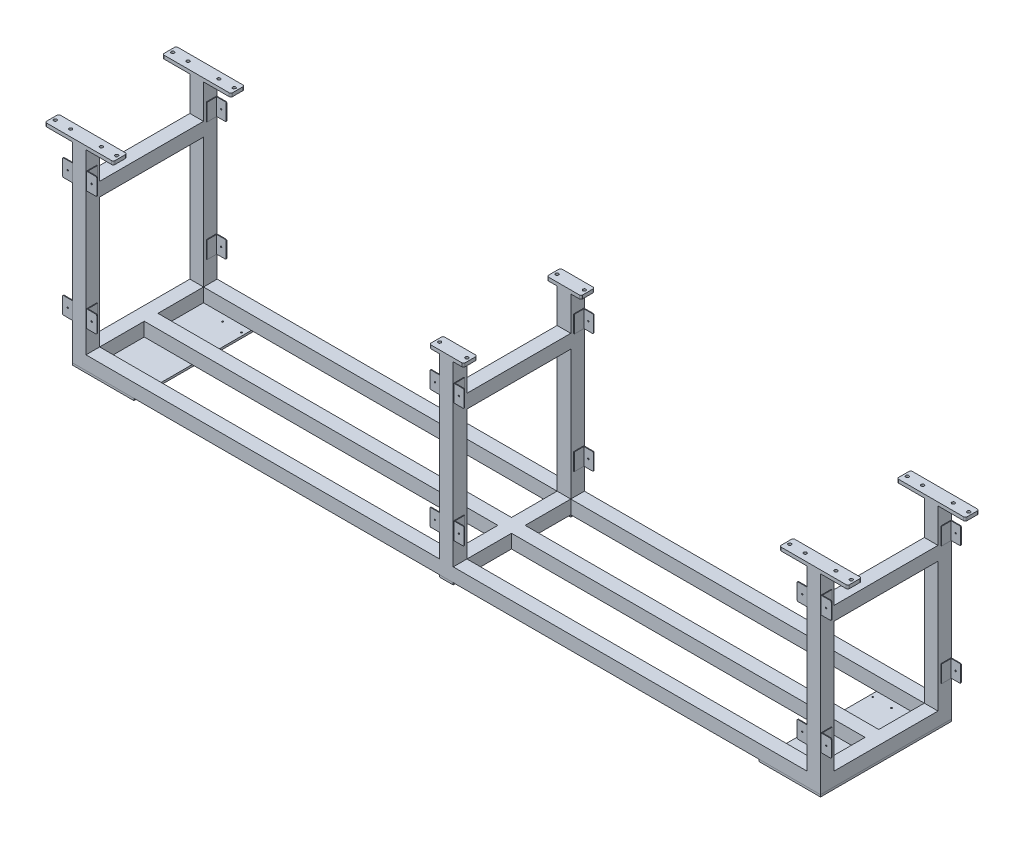
SolidWorks part; units mm, degrees
ref_plane "前视基准面" through (0, 0, 0) normal (0, 0, 1) x (1, 0, 0)
ref_plane "上视基准面" through (0, 0, 0) normal (0, 1, 0) x (1, 0, 0)
ref_plane "右视基准面" through (0, 0, 0) normal (1, 0, 0) x (0, 0, -1)
sketch "草图1" plane through (0, 0, 0) normal (0, 0, 1) x (1, 0, 0)
  line L0 (-81.7263, -196.6753) -> (953.2737, -196.6753)
  line L1 (-81.7263, -156.6753) -> (953.2737, -156.6753)
  line L2 (-81.7263, -161.6753) -> (953.2737, -161.6753) construction
  line L3 (-81.7263, -191.6753) -> (953.2737, -191.6753) construction
  line L4 (-121.7263, -196.6753) -> (-1186.7263, -196.6753)
  line L5 (-121.7263, -156.6753) -> (-1186.7263, -156.6753)
  line L6 (-121.7263, -161.6753) -> (-1186.7263, -161.6753) construction
  line L7 (-121.7263, -191.6753) -> (-1186.7263, -191.6753) construction
  line L8 (-1186.7263, -196.6753) -> (-1196.7263, -196.6753)
  line L9 (-1196.7263, -196.6753) -> (-1196.7263, -156.6753)
  line L10 (-1186.7263, -156.6753) -> (-1196.7263, -156.6753)
  line L11 (993.2737, -196.6753) -> (953.2737, -196.6753)
  line L12 (973.2737, -176.2036) -> (973.2737, -230.0906) construction
  line L13 (993.2737, -196.6753) -> (813.2737, -196.6753)
  line L14 (813.2737, -196.6753) -> (813.2737, -202.6753)
  line L15 (813.2737, -202.6753) -> (993.2737, -202.6753)
  line L16 (993.2737, -196.6753) -> (993.2737, -202.6753)
  line L17 (966.3455, -204.6753) -> (966.3455, -216.6753)
  line L18 (980.2019, -204.6753) -> (980.2019, -216.6753)
  line L19 (962.8814, -218.6753) -> (983.666, -218.6753)
  line L20 (959.4173, -204.6753) -> (959.4173, -216.6753)
  line L21 (987.1301, -204.6753) -> (987.1301, -216.6753)
  line L22 (962.8814, -202.6753) -> (983.666, -202.6753)
  line L23 (-1196.7263, -196.6753) -> (-1156.7263, -196.6753)
  line L24 (-1196.7263, -196.6753) -> (-1016.7263, -196.6753)
  line L25 (-1016.7263, -196.6753) -> (-1016.7263, -202.6753)
  line L26 (-1016.7263, -202.6753) -> (-1196.7263, -202.6753)
  line L27 (-1196.7263, -196.6753) -> (-1196.7263, -202.6753)
  line L28 (-1169.7981, -204.6753) -> (-1169.7981, -216.6753)
  line L29 (-1183.6545, -204.6753) -> (-1183.6545, -216.6753)
  line L30 (-1166.334, -218.6753) -> (-1187.1186, -218.6753)
  line L31 (-1162.8699, -204.6753) -> (-1162.8699, -216.6753)
  line L32 (-1190.5827, -204.6753) -> (-1190.5827, -216.6753)
  line L33 (-1166.334, -202.6753) -> (-1187.1186, -202.6753)
  line L34 (-1146.5223, -176.6753) -> (-1216.0939, -176.6753) construction
  line L35 (943.0697, -176.6753) -> (1012.6413, -176.6753) construction
  spline S0 degree 3 poles (959.4173, -216.6753) (960.572, -217.6753) (962.8814, -219.6753) (965.1908, -217.6753) (966.3455, -216.6753) knots 0 0 0 0 0.5 1 1 1 1
  spline S1 degree 3 poles (966.3455, -216.6753) (968.6549, -217.6753) (973.2737, -219.6753) (977.8925, -217.6753) (980.2019, -216.6753) knots 0 0 0 0 0.5 1 1 1 1
  spline S2 degree 3 poles (987.1301, -216.6753) (985.9754, -217.6753) (983.666, -219.6753) (981.3566, -217.6753) (980.2019, -216.6753) knots 0 0 0 0 0.5 1 1 1 1
  spline S3 degree 3 poles (966.3455, -204.6753) (968.6549, -203.6753) (973.2737, -201.6753) (977.8925, -203.6753) (980.2019, -204.6753) knots 0 0 0 0 0.5 1 1 1 1
  spline S4 degree 3 poles (959.4173, -204.6753) (960.572, -203.6753) (962.8814, -201.6753) (965.1908, -203.6753) (966.3455, -204.6753) knots 0 0 0 0 0.5 1 1 1 1
  spline S5 degree 3 poles (987.1301, -204.6753) (985.9754, -203.6753) (983.666, -201.6753) (981.3566, -203.6753) (980.2019, -204.6753) knots 0 0 0 0 0.5 1 1 1 1
  spline S6 degree 3 poles (-1162.8699, -216.6753) (-1164.0246, -217.6753) (-1166.334, -219.6753) (-1168.6434, -217.6753) (-1169.7981, -216.6753) knots 0 0 0 0 0.5 1 1 1 1
  spline S7 degree 3 poles (-1169.7981, -216.6753) (-1172.1075, -217.6753) (-1176.7263, -219.6753) (-1181.3451, -217.6753) (-1183.6545, -216.6753) knots 0 0 0 0 0.5 1 1 1 1
  spline S8 degree 3 poles (-1190.5827, -216.6753) (-1189.428, -217.6753) (-1187.1186, -219.6753) (-1184.8092, -217.6753) (-1183.6545, -216.6753) knots 0 0 0 0 0.5 1 1 1 1
  spline S9 degree 3 poles (-1169.7981, -204.6753) (-1172.1075, -203.6753) (-1176.7263, -201.6753) (-1181.3451, -203.6753) (-1183.6545, -204.6753) knots 0 0 0 0 0.5 1 1 1 1
  spline S10 degree 3 poles (-1162.8699, -204.6753) (-1164.0246, -203.6753) (-1166.334, -201.6753) (-1168.6434, -203.6753) (-1169.7981, -204.6753) knots 0 0 0 0 0.5 1 1 1 1
  spline S11 degree 3 poles (-1190.5827, -204.6753) (-1189.428, -203.6753) (-1187.1186, -201.6753) (-1184.8092, -203.6753) (-1183.6545, -204.6753) knots 0 0 0 0 0.5 1 1 1 1
  line B0 (-121.7263, 363.3247) -> (-121.7263, -196.6753)
  line B1 (-116.7263, 363.3247) -> (-116.7263, -196.6753) construction
  line B2 (-121.7263, -196.6753) -> (-81.7263, -196.6753)
  line B3 (-116.7263, -186.6753) -> (-86.7263, -186.6753) construction
  line B4 (-81.7263, -196.6753) -> (-81.7263, 363.3247)
  line B5 (-86.7263, -196.6753) -> (-86.7263, 363.3247) construction
  line B6 (-151.7263, 373.3247) -> (-51.7263, 373.3247)
  line B7 (-151.7263, 363.3247) -> (-51.7263, 363.3247)
  line B8 (-151.7263, 373.3247) -> (-151.7263, 363.3247)
  line B9 (-51.7263, 373.3247) -> (-51.7263, 363.3247)
  line B10 (-101.7263, -176.2036) -> (-101.7263, -206.1494) construction
  line B11 (-109.7263, -186.6753) -> (-109.7263, -196.6753) construction
  line B12 (-108.2263, -186.6753) -> (-108.2263, -196.6753) construction
  line B13 (-93.7263, -186.6753) -> (-93.7263, -196.6753) construction
  line B14 (-95.2263, -186.6753) -> (-95.2263, -196.6753) construction
  line B15 (-61.7263, 352.831) -> (-61.7263, 383.9585) construction
  line B16 (-141.7263, 352.831) -> (-141.7263, 383.9585) construction
  line B17 (-121.7263, -156.6753) -> (-81.7263, -156.6753) construction
  line B18 (-81.7263, -156.6753) -> (-81.7263, -196.6753) construction
  line B19 (-81.7263, -196.6753) -> (-121.7263, -196.6753) construction
  line B20 (-121.7263, -196.6753) -> (-121.7263, -156.6753) construction
  line B21 (-116.7263, -161.6753) -> (-86.7263, -161.6753) construction
  line B22 (-86.7263, -161.6753) -> (-86.7263, -191.6753) construction
  line B23 (-86.7263, -191.6753) -> (-116.7263, -191.6753) construction
  line B24 (-116.7263, -191.6753) -> (-116.7263, -161.6753) construction
  line B25 (-121.7263, 263.3247) -> (-81.7263, 263.3247) construction
  line B26 (-81.7263, 263.3247) -> (-81.7263, 223.3247) construction
  line B27 (-81.7263, 223.3247) -> (-121.7263, 223.3247) construction
  line B28 (-121.7263, 223.3247) -> (-121.7263, 263.3247) construction
  line B29 (-116.7263, 258.3247) -> (-86.7263, 258.3247) construction
  line B30 (-86.7263, 258.3247) -> (-86.7263, 228.3247) construction
  line B31 (-86.7263, 228.3247) -> (-116.7263, 228.3247) construction
  line B32 (-116.7263, 228.3247) -> (-116.7263, 258.3247) construction
  line B33 (-108.7263, -196.6753) -> (-108.7263, -268.6753)
  line B34 (-109.7263, -196.6753) -> (-109.7263, -268.6753)
  line B35 (-94.7263, -196.6753) -> (-94.7263, -268.6753)
  line B36 (-93.7263, -196.6753) -> (-93.7263, -268.6753)
  line B37 (-131.7263, -287.6753) -> (-131.7263, -288.6753)
  line B38 (-71.7263, -287.6753) -> (-71.7263, -288.6753)
  line B39 (-71.7263, -288.6753) -> (-131.7263, -288.6753)
  line B40 (-71.7263, -287.6753) -> (-131.7263, -287.6753)
  line B41 (-84.7263, -278.6753) -> (-118.7263, -278.6753)
  line B42 (-114.7263, -270.1755) -> (-114.7263, -277.1751)
  line B43 (-109.2263, -270.1753) -> (-109.2263, -277.1755)
  line B44 (-91.3223, -268.6753) -> (-111.944, -268.6753)
  line B45 (-91.4763, -268.6753) -> (-111.9762, -268.6753)
  line B46 (-94.2263, -270.1753) -> (-94.2263, -277.1753)
  line B47 (-88.7263, -270.1753) -> (-88.7263, -277.1753)
  line B48 (-109.7263, -196.6753) -> (-93.7263, -196.6753)
  arc B49 (-94.2263, -277.1753) -> (-88.7263, -277.1753) centre (-91.4763, -275.4045) ccw
  arc B50 (-76.7263, -287.6753) -> (-84.7263, -278.6753) centre (-95.3954, -296.2145) ccw
  arc B51 (-109.2263, -277.1753) -> (-94.2263, -277.1753) centre (-101.7263, -259.1753) ccw
  arc B52 (-114.7262, -277.1753) -> (-109.2262, -277.1753) centre (-111.9762, -275.4045) ccw
  arc B53 (-118.7261, -278.6753) -> (-126.7261, -287.6753) centre (-108.0569, -296.2145) ccw
  arc B54 (-109.2262, -270.1753) -> (-114.7262, -270.1753) centre (-111.9762, -271.9461) ccw
  arc B55 (-94.2263, -270.1753) -> (-109.2263, -270.1753) centre (-101.7263, -288.1753) ccw
  arc B56 (-88.7263, -270.1753) -> (-94.2263, -270.1753) centre (-91.4763, -271.9461) ccw
  line B57 (980.2737, -218.6753) -> (980.2737, -268.6753)
  line B58 (981.2737, -218.6753) -> (981.2737, -268.6753)
  line B59 (966.2737, -218.6753) -> (966.2737, -268.6753)
  line B60 (965.2737, -218.6753) -> (965.2737, -268.6753)
  line B61 (1003.2737, -287.6753) -> (1003.2737, -288.6753)
  line B62 (943.2737, -287.6753) -> (943.2737, -288.6753)
  line B63 (943.2737, -288.6753) -> (1003.2737, -288.6753)
  line B64 (943.2737, -287.6753) -> (1003.2737, -287.6753)
  line B65 (956.2737, -278.6753) -> (990.2737, -278.6753)
  line B66 (986.2737, -270.1755) -> (986.2737, -277.1751)
  line B67 (980.7737, -270.1753) -> (980.7737, -277.1755)
  line B68 (962.8697, -268.6753) -> (983.4914, -268.6753)
  line B69 (963.0237, -268.6753) -> (983.5236, -268.6753)
  line B70 (965.7737, -270.1753) -> (965.7737, -277.1753)
  line B71 (960.2737, -270.1753) -> (960.2737, -277.1753)
  line B72 (981.2737, -218.6753) -> (965.2737, -218.6753)
  arc B73 (960.2737, -277.1753) -> (965.7737, -277.1753) centre (963.0237, -275.4045) ccw
  arc B74 (956.2737, -278.6753) -> (948.2737, -287.6753) centre (966.9428, -296.2145) ccw
  arc B75 (965.7737, -277.1753) -> (980.7737, -277.1753) centre (973.2737, -259.1753) ccw
  arc B76 (980.7736, -277.1753) -> (986.2736, -277.1753) centre (983.5236, -275.4045) ccw
  arc B77 (998.2735, -287.6753) -> (990.2735, -278.6753) centre (979.6044, -296.2145) ccw
  arc B78 (986.2736, -270.1753) -> (980.7736, -270.1753) centre (983.5236, -271.9461) ccw
  arc B79 (980.7737, -270.1753) -> (965.7737, -270.1753) centre (973.2737, -288.1753) ccw
  arc B80 (965.7737, -270.1753) -> (960.2737, -270.1753) centre (963.0237, -271.9461) ccw
  line B81 (893.2737, -229.6753) -> (893.2737, -223.6753)
  line B82 (888.2737, -218.6753) -> (838.2737, -218.6753)
  line B83 (828.3708, -223.6753) -> (827.5097, -229.6753)
  line B84 (903.2737, -208.6753) -> (813.2737, -208.6753)
  line B85 (813.2737, -208.6753) -> (813.2737, -202.6753)
  line B86 (813.2737, -202.6753) -> (903.2737, -202.6753)
  line B87 (903.2737, -202.6753) -> (903.2737, -208.6753)
  line B88 (888.2737, -208.6753) -> (888.2737, -218.6753)
  line B89 (888.2737, -218.6753) -> (838.2737, -218.6753)
  line B90 (838.2737, -218.6753) -> (838.2737, -208.6753)
  line B91 (838.2737, -208.6753) -> (888.2737, -208.6753)
  line B92 (893.2737, -229.6753) -> (893.2737, -223.6753)
  line B93 (888.2737, -218.6753) -> (838.2737, -218.6753)
  line B94 (828.3708, -223.6753) -> (827.5097, -229.6753)
  line B95 (903.2737, -208.6753) -> (813.2737, -208.6753)
  line B96 (813.2737, -208.6753) -> (813.2737, -202.6753)
  line B97 (813.2737, -202.6753) -> (903.2737, -202.6753)
  line B98 (903.2737, -202.6753) -> (903.2737, -208.6753)
  line B99 (888.2737, -208.6753) -> (888.2737, -218.6753)
  line B100 (888.2737, -218.6753) -> (838.2737, -218.6753)
  line B101 (838.2737, -218.6753) -> (838.2737, -208.6753)
  line B102 (838.2737, -208.6753) -> (888.2737, -208.6753)
  arc B103 (893.2737, -223.6753) -> (888.2737, -218.6753) centre (888.2737, -223.6753) ccw
  arc B104 (838.2737, -218.6753) -> (828.3708, -223.6753) centre (837.7267, -229.8987) ccw
  arc B105 (826.9708, -240.4435) -> (859.8834, -242.2847) centre (842.7943, -252.6753) ccw
  arc B106 (827.9504, -226.6051) -> (866.767, -234.6389) centre (842.7943, -252.6753) ccw
  circle B107 centre (842.7943, -252.6753) radius 6
  arc B108 (893.2737, -223.6753) -> (888.2737, -218.6753) centre (888.2737, -223.6753) ccw
  arc B109 (838.2737, -218.6753) -> (828.3708, -223.6753) centre (837.7267, -229.8987) ccw
  arc B110 (826.9708, -240.4435) -> (859.8834, -242.2847) centre (842.7943, -252.6753) ccw
  arc B111 (827.9504, -226.6051) -> (866.767, -234.6389) centre (842.7943, -252.6753) ccw
  circle B112 centre (842.7943, -252.6753) radius 6
  spline B113 degree 3 poles (893.2737, -229.6753) (889.5179, -229.4713) (877.6067, -228.8243) (856.7832, -237.1379) (858.2534, -263.4691) (830.1026, -264.2073) (826.3694, -244.5927) (827.1435, -234.466) (827.5097, -229.6753) knots 0 0 0 0 0.107435 0.340721 0.514208 0.707478 0.861613 1 1 1 1
  spline B114 degree 3 poles (893.2737, -229.6753) (889.5179, -229.4713) (877.6067, -228.8243) (856.7832, -237.1379) (858.2534, -263.4691) (830.1026, -264.2073) (826.3694, -244.5927) (827.1435, -234.466) (827.5097, -229.6753) knots 0 0 0 0 0.107435 0.340721 0.514208 0.707478 0.861613 1 1 1 1
  line B115 (-81.7263, 308.3247) -> (-54.7263, 308.3247)
  line B116 (-51.7263, 305.3247) -> (-51.7263, 261.3247)
  line B117 (-54.7263, 258.3247) -> (-81.7263, 258.3247)
  line B118 (-81.7263, 258.3247) -> (-81.7263, 308.3247)
  line B119 (-79.7263, 258.3247) -> (-79.7263, 308.3247) construction
  arc B120 (-51.7263, 305.3247) -> (-54.7263, 308.3247) centre (-54.7263, 305.3247) ccw
  arc B121 (-54.7263, 258.3247) -> (-51.7263, 261.3247) centre (-54.7263, 261.3247) ccw
  arc B122 (-64.2263, 283.3247) -> (-66.7263, 280.8247) centre (-66.7263, 283.3247) ccw
  circle B123 centre (-66.7263, 283.3247) radius 2
  line B124 (-81.7263, -40.6753) -> (-54.7263, -40.6753)
  line B125 (-51.7263, -43.6753) -> (-51.7263, -87.6753)
  line B126 (-54.7263, -90.6753) -> (-81.7263, -90.6753)
  line B127 (-81.7263, -90.6753) -> (-81.7263, -40.6753)
  line B128 (-79.7263, -90.6753) -> (-79.7263, -40.6753) construction
  arc B129 (-51.7263, -43.6753) -> (-54.7263, -40.6753) centre (-54.7263, -43.6753) ccw
  arc B130 (-54.7263, -90.6753) -> (-51.7263, -87.6753) centre (-54.7263, -87.6753) ccw
  arc B131 (-64.2263, -65.6753) -> (-66.7263, -68.1753) centre (-66.7263, -65.6753) ccw
  circle B132 centre (-66.7263, -65.6753) radius 2
  line B133 (-121.7263, 308.3247) -> (-148.7263, 308.3247)
  line B134 (-151.7263, 305.3247) -> (-151.7263, 261.3247)
  line B135 (-148.7263, 258.3247) -> (-121.7263, 258.3247)
  line B136 (-121.7263, 258.3247) -> (-121.7263, 308.3247)
  line B137 (-123.7263, 258.3247) -> (-123.7263, 308.3247) construction
  arc B138 (-148.7263, 308.3247) -> (-151.7263, 305.3247) centre (-148.7263, 305.3247) ccw
  arc B139 (-151.7263, 261.3247) -> (-148.7263, 258.3247) centre (-148.7263, 261.3247) ccw
  arc B140 (-136.7263, 280.8247) -> (-139.2263, 283.3247) centre (-136.7263, 283.3247) ccw
  circle B141 centre (-136.7263, 283.3247) radius 2
  line B142 (-121.7263, -40.6753) -> (-148.7263, -40.6753)
  line B143 (-151.7263, -43.6753) -> (-151.7263, -87.6753)
  line B144 (-148.7263, -90.6753) -> (-121.7263, -90.6753)
  line B145 (-121.7263, -90.6753) -> (-121.7263, -40.6753)
  line B146 (-123.7263, -90.6753) -> (-123.7263, -40.6753) construction
  arc B147 (-148.7263, -40.6753) -> (-151.7263, -43.6753) centre (-148.7263, -43.6753) ccw
  arc B148 (-151.7263, -87.6753) -> (-148.7263, -90.6753) centre (-148.7263, -87.6753) ccw
  arc B149 (-136.7263, -68.1753) -> (-139.2263, -65.6753) centre (-136.7263, -65.6753) ccw
  circle B150 centre (-136.7263, -65.6753) radius 2
  line B151 (953.2737, 363.3247) -> (953.2737, -196.6753)
  line B152 (958.2737, 363.3247) -> (958.2737, -196.6753) construction
  line B153 (953.2737, -196.6753) -> (993.2737, -196.6753)
  line B154 (958.2737, -186.6753) -> (988.2737, -186.6753) construction
  line B155 (993.2737, -196.6753) -> (993.2737, 363.3247)
  line B156 (988.2737, -196.6753) -> (988.2737, 363.3247) construction
  line B157 (873.2737, 373.3247) -> (1073.2737, 373.3247)
  line B158 (873.2737, 363.3247) -> (1073.2737, 363.3247)
  line B159 (873.2737, 373.3247) -> (873.2737, 363.3247)
  line B160 (1073.2737, 373.3247) -> (1073.2737, 363.3247)
  line B161 (973.2737, -176.2036) -> (973.2737, -206.1494) construction
  line B162 (965.2737, -186.6753) -> (965.2737, -196.6753) construction
  line B163 (966.7737, -186.6753) -> (966.7737, -196.6753) construction
  line B164 (981.2737, -186.6753) -> (981.2737, -196.6753) construction
  line B165 (979.7737, -186.6753) -> (979.7737, -196.6753) construction
  line B166 (1063.2737, 352.831) -> (1063.2737, 383.9585) construction
  line B167 (883.2737, 352.831) -> (883.2737, 383.9585) construction
  line B168 (1018.2737, 352.831) -> (1018.2737, 383.9585) construction
  line B169 (928.2737, 352.831) -> (928.2737, 383.9585) construction
  line B170 (953.2737, 263.3247) -> (993.2737, 263.3247) construction
  line B171 (993.2737, 263.3247) -> (993.2737, 223.3247) construction
  line B172 (993.2737, 223.3247) -> (953.2737, 223.3247) construction
  line B173 (953.2737, 223.3247) -> (953.2737, 263.3247) construction
  line B174 (958.2737, 258.3247) -> (988.2737, 258.3247) construction
  line B175 (988.2737, 258.3247) -> (988.2737, 228.3247) construction
  line B176 (988.2737, 228.3247) -> (958.2737, 228.3247) construction
  line B177 (958.2737, 228.3247) -> (958.2737, 258.3247) construction
  line B178 (953.2737, -156.6753) -> (993.2737, -156.6753) construction
  line B179 (993.2737, -156.6753) -> (993.2737, -196.6753) construction
  line B180 (993.2737, -196.6753) -> (953.2737, -196.6753) construction
  line B181 (953.2737, -196.6753) -> (953.2737, -156.6753) construction
  line B182 (958.2737, -161.6753) -> (988.2737, -161.6753) construction
  line B183 (988.2737, -161.6753) -> (988.2737, -191.6753) construction
  line B184 (988.2737, -191.6753) -> (958.2737, -191.6753) construction
  line B185 (958.2737, -191.6753) -> (958.2737, -161.6753) construction
  line B186 (993.2737, 308.3247) -> (1020.2737, 308.3247)
  line B187 (1023.2737, 305.3247) -> (1023.2737, 261.3247)
  line B188 (1020.2737, 258.3247) -> (993.2737, 258.3247)
  line B189 (993.2737, 258.3247) -> (993.2737, 308.3247)
  line B190 (995.2737, 258.3247) -> (995.2737, 308.3247) construction
  arc B191 (1023.2737, 305.3247) -> (1020.2737, 308.3247) centre (1020.2737, 305.3247) ccw
  arc B192 (1020.2737, 258.3247) -> (1023.2737, 261.3247) centre (1020.2737, 261.3247) ccw
  arc B193 (1010.7737, 283.3247) -> (1008.2737, 280.8247) centre (1008.2737, 283.3247) ccw
  circle B194 centre (1008.2737, 283.3247) radius 2
  line B195 (993.2737, -40.6753) -> (1020.2737, -40.6753)
  line B196 (1023.2737, -43.6753) -> (1023.2737, -87.6753)
  line B197 (1020.2737, -90.6753) -> (993.2737, -90.6753)
  line B198 (993.2737, -90.6753) -> (993.2737, -40.6753)
  line B199 (995.2737, -90.6753) -> (995.2737, -40.6753) construction
  arc B200 (1023.2737, -43.6753) -> (1020.2737, -40.6753) centre (1020.2737, -43.6753) ccw
  arc B201 (1020.2737, -90.6753) -> (1023.2737, -87.6753) centre (1020.2737, -87.6753) ccw
  arc B202 (1010.7737, -65.6753) -> (1008.2737, -68.1753) centre (1008.2737, -65.6753) ccw
  circle B203 centre (1008.2737, -65.6753) radius 2
  line B204 (953.2737, 308.3247) -> (926.2737, 308.3247)
  line B205 (923.2737, 305.3247) -> (923.2737, 261.3247)
  line B206 (926.2737, 258.3247) -> (953.2737, 258.3247)
  line B207 (953.2737, 258.3247) -> (953.2737, 308.3247)
  line B208 (951.2737, 258.3247) -> (951.2737, 308.3247) construction
  arc B209 (926.2737, 308.3247) -> (923.2737, 305.3247) centre (926.2737, 305.3247) ccw
  arc B210 (923.2737, 261.3247) -> (926.2737, 258.3247) centre (926.2737, 261.3247) ccw
  arc B211 (938.2737, 280.8247) -> (935.7737, 283.3247) centre (938.2737, 283.3247) ccw
  circle B212 centre (938.2737, 283.3247) radius 2
  line B213 (953.2737, -40.6753) -> (926.2737, -40.6753)
  line B214 (923.2737, -43.6753) -> (923.2737, -87.6753)
  line B215 (926.2737, -90.6753) -> (953.2737, -90.6753)
  line B216 (953.2737, -90.6753) -> (953.2737, -40.6753)
  line B217 (951.2737, -90.6753) -> (951.2737, -40.6753) construction
  arc B218 (926.2737, -40.6753) -> (923.2737, -43.6753) centre (926.2737, -43.6753) ccw
  arc B219 (923.2737, -87.6753) -> (926.2737, -90.6753) centre (926.2737, -87.6753) ccw
  arc B220 (938.2737, -68.1753) -> (935.7737, -65.6753) centre (938.2737, -65.6753) ccw
  circle B221 centre (938.2737, -65.6753) radius 2
  line B222 (-1183.7263, -218.6753) -> (-1183.7263, -268.6753)
  line B223 (-1184.7263, -218.6753) -> (-1184.7263, -268.6753)
  line B224 (-1169.7263, -218.6753) -> (-1169.7263, -268.6753)
  line B225 (-1168.7263, -218.6753) -> (-1168.7263, -268.6753)
  line B226 (-1206.7263, -287.6753) -> (-1206.7263, -288.6753)
  line B227 (-1146.7263, -287.6753) -> (-1146.7263, -288.6753)
  line B228 (-1146.7263, -288.6753) -> (-1206.7263, -288.6753)
  line B229 (-1146.7263, -287.6753) -> (-1206.7263, -287.6753)
  line B230 (-1159.7263, -278.6753) -> (-1193.7263, -278.6753)
  line B231 (-1189.7263, -270.1755) -> (-1189.7263, -277.1751)
  line B232 (-1184.2263, -270.1753) -> (-1184.2263, -277.1755)
  line B233 (-1166.3223, -268.6753) -> (-1186.944, -268.6753)
  line B234 (-1166.4763, -268.6753) -> (-1186.9762, -268.6753)
  line B235 (-1169.2263, -270.1753) -> (-1169.2263, -277.1753)
  line B236 (-1163.7263, -270.1753) -> (-1163.7263, -277.1753)
  line B237 (-1184.7263, -218.6753) -> (-1168.7263, -218.6753)
  arc B238 (-1169.2263, -277.1753) -> (-1163.7263, -277.1753) centre (-1166.4763, -275.4045) ccw
  arc B239 (-1151.7263, -287.6753) -> (-1159.7263, -278.6753) centre (-1170.3954, -296.2145) ccw
  arc B240 (-1184.2263, -277.1753) -> (-1169.2263, -277.1753) centre (-1176.7263, -259.1753) ccw
  arc B241 (-1189.7262, -277.1753) -> (-1184.2262, -277.1753) centre (-1186.9762, -275.4045) ccw
  arc B242 (-1193.7261, -278.6753) -> (-1201.7261, -287.6753) centre (-1183.0569, -296.2145) ccw
  arc B243 (-1184.2262, -270.1753) -> (-1189.7262, -270.1753) centre (-1186.9762, -271.9461) ccw
  arc B244 (-1169.2263, -270.1753) -> (-1184.2263, -270.1753) centre (-1176.7263, -288.1753) ccw
  arc B245 (-1163.7263, -270.1753) -> (-1169.2263, -270.1753) centre (-1166.4763, -271.9461) ccw
  line B246 (-1096.7263, -229.6753) -> (-1096.7263, -223.6753)
  line B247 (-1091.7263, -218.6753) -> (-1041.7263, -218.6753)
  line B248 (-1031.8234, -223.6753) -> (-1030.9623, -229.6753)
  line B249 (-1106.7263, -208.6753) -> (-1016.7263, -208.6753)
  line B250 (-1016.7263, -208.6753) -> (-1016.7263, -202.6753)
  line B251 (-1016.7263, -202.6753) -> (-1106.7263, -202.6753)
  line B252 (-1106.7263, -202.6753) -> (-1106.7263, -208.6753)
  line B253 (-1091.7263, -208.6753) -> (-1091.7263, -218.6753)
  line B254 (-1091.7263, -218.6753) -> (-1041.7263, -218.6753)
  line B255 (-1041.7263, -218.6753) -> (-1041.7263, -208.6753)
  line B256 (-1041.7263, -208.6753) -> (-1091.7263, -208.6753)
  line B257 (-1096.7263, -229.6753) -> (-1096.7263, -223.6753)
  line B258 (-1091.7263, -218.6753) -> (-1041.7263, -218.6753)
  line B259 (-1031.8234, -223.6753) -> (-1030.9623, -229.6753)
  line B260 (-1106.7263, -208.6753) -> (-1016.7263, -208.6753)
  line B261 (-1016.7263, -208.6753) -> (-1016.7263, -202.6753)
  line B262 (-1016.7263, -202.6753) -> (-1106.7263, -202.6753)
  line B263 (-1106.7263, -202.6753) -> (-1106.7263, -208.6753)
  line B264 (-1091.7263, -208.6753) -> (-1091.7263, -218.6753)
  line B265 (-1091.7263, -218.6753) -> (-1041.7263, -218.6753)
  line B266 (-1041.7263, -218.6753) -> (-1041.7263, -208.6753)
  line B267 (-1041.7263, -208.6753) -> (-1091.7263, -208.6753)
  arc B268 (-1091.7263, -218.6753) -> (-1096.7263, -223.6753) centre (-1091.7263, -223.6753) ccw
  arc B269 (-1031.8234, -223.6753) -> (-1041.7263, -218.6753) centre (-1041.1793, -229.8987) ccw
  arc B270 (-1063.336, -242.2847) -> (-1030.4234, -240.4435) centre (-1046.2469, -252.6753) ccw
  arc B271 (-1070.2196, -234.6389) -> (-1031.4029, -226.6051) centre (-1046.2469, -252.6753) ccw
  circle B272 centre (-1046.2469, -252.6753) radius 6
  arc B273 (-1091.7263, -218.6753) -> (-1096.7263, -223.6753) centre (-1091.7263, -223.6753) ccw
  arc B274 (-1031.8234, -223.6753) -> (-1041.7263, -218.6753) centre (-1041.1793, -229.8987) ccw
  arc B275 (-1063.336, -242.2847) -> (-1030.4234, -240.4435) centre (-1046.2469, -252.6753) ccw
  arc B276 (-1070.2196, -234.6389) -> (-1031.4029, -226.6051) centre (-1046.2469, -252.6753) ccw
  circle B277 centre (-1046.2469, -252.6753) radius 6
  spline B278 degree 3 poles (-1096.7263, -229.6753) (-1092.9705, -229.4713) (-1081.0593, -228.8243) (-1060.2358, -237.1379) (-1061.7059, -263.4691) (-1033.5552, -264.2073) (-1029.822, -244.5927) (-1030.5961, -234.466) (-1030.9623, -229.6753) knots 0 0 0 0 0.107435 0.340721 0.514208 0.707478 0.861613 1 1 1 1
  spline B279 degree 3 poles (-1096.7263, -229.6753) (-1092.9705, -229.4713) (-1081.0593, -228.8243) (-1060.2358, -237.1379) (-1061.7059, -263.4691) (-1033.5552, -264.2073) (-1029.822, -244.5927) (-1030.5961, -234.466) (-1030.9623, -229.6753) knots 0 0 0 0 0.107435 0.340721 0.514208 0.707478 0.861613 1 1 1 1
  line B280 (-1156.7263, 363.3247) -> (-1156.7263, -196.6753)
  line B281 (-1161.7263, 363.3247) -> (-1161.7263, -196.6753) construction
  line B282 (-1156.7263, -196.6753) -> (-1196.7263, -196.6753)
  line B283 (-1161.7263, -186.6753) -> (-1191.7263, -186.6753) construction
  line B284 (-1196.7263, -196.6753) -> (-1196.7263, 363.3247)
  line B285 (-1191.7263, -196.6753) -> (-1191.7263, 363.3247) construction
  line B286 (-1076.7263, 373.3247) -> (-1276.7263, 373.3247)
  line B287 (-1076.7263, 363.3247) -> (-1276.7263, 363.3247)
  line B288 (-1076.7263, 373.3247) -> (-1076.7263, 363.3247)
  line B289 (-1276.7263, 373.3247) -> (-1276.7263, 363.3247)
  line B290 (-1176.7263, -176.2036) -> (-1176.7263, -206.1494) construction
  line B291 (-1168.7263, -186.6753) -> (-1168.7263, -196.6753) construction
  line B292 (-1170.2263, -186.6753) -> (-1170.2263, -196.6753) construction
  line B293 (-1184.7263, -186.6753) -> (-1184.7263, -196.6753) construction
  line B294 (-1183.2263, -186.6753) -> (-1183.2263, -196.6753) construction
  line B295 (-1266.7263, 352.831) -> (-1266.7263, 383.9585) construction
  line B296 (-1086.7263, 352.831) -> (-1086.7263, 383.9585) construction
  line B297 (-1221.7263, 352.831) -> (-1221.7263, 383.9585) construction
  line B298 (-1131.7263, 352.831) -> (-1131.7263, 383.9585) construction
  line B299 (-1156.7263, 263.3247) -> (-1196.7263, 263.3247) construction
  line B300 (-1196.7263, 263.3247) -> (-1196.7263, 223.3247) construction
  line B301 (-1196.7263, 223.3247) -> (-1156.7263, 223.3247) construction
  line B302 (-1156.7263, 223.3247) -> (-1156.7263, 263.3247) construction
  line B303 (-1161.7263, 258.3247) -> (-1191.7263, 258.3247) construction
  line B304 (-1191.7263, 258.3247) -> (-1191.7263, 228.3247) construction
  line B305 (-1191.7263, 228.3247) -> (-1161.7263, 228.3247) construction
  line B306 (-1161.7263, 228.3247) -> (-1161.7263, 258.3247) construction
  line B307 (-1156.7263, -156.6753) -> (-1196.7263, -156.6753) construction
  line B308 (-1196.7263, -156.6753) -> (-1196.7263, -196.6753) construction
  line B309 (-1196.7263, -196.6753) -> (-1156.7263, -196.6753) construction
  line B310 (-1156.7263, -196.6753) -> (-1156.7263, -156.6753) construction
  line B311 (-1161.7263, -161.6753) -> (-1191.7263, -161.6753) construction
  line B312 (-1191.7263, -161.6753) -> (-1191.7263, -191.6753) construction
  line B313 (-1191.7263, -191.6753) -> (-1161.7263, -191.6753) construction
  line B314 (-1161.7263, -191.6753) -> (-1161.7263, -161.6753) construction
  line B315 (-1196.7263, 308.3247) -> (-1223.7263, 308.3247)
  line B316 (-1226.7263, 305.3247) -> (-1226.7263, 261.3247)
  line B317 (-1223.7263, 258.3247) -> (-1196.7263, 258.3247)
  line B318 (-1196.7263, 258.3247) -> (-1196.7263, 308.3247)
  line B319 (-1198.7263, 258.3247) -> (-1198.7263, 308.3247) construction
  arc B320 (-1223.7263, 308.3247) -> (-1226.7263, 305.3247) centre (-1223.7263, 305.3247) ccw
  arc B321 (-1226.7263, 261.3247) -> (-1223.7263, 258.3247) centre (-1223.7263, 261.3247) ccw
  arc B322 (-1211.7263, 280.8247) -> (-1214.2263, 283.3247) centre (-1211.7263, 283.3247) ccw
  circle B323 centre (-1211.7263, 283.3247) radius 2
  line B324 (-1196.7263, -40.6753) -> (-1223.7263, -40.6753)
  line B325 (-1226.7263, -43.6753) -> (-1226.7263, -87.6753)
  line B326 (-1223.7263, -90.6753) -> (-1196.7263, -90.6753)
  line B327 (-1196.7263, -90.6753) -> (-1196.7263, -40.6753)
  line B328 (-1198.7263, -90.6753) -> (-1198.7263, -40.6753) construction
  arc B329 (-1223.7263, -40.6753) -> (-1226.7263, -43.6753) centre (-1223.7263, -43.6753) ccw
  arc B330 (-1226.7263, -87.6753) -> (-1223.7263, -90.6753) centre (-1223.7263, -87.6753) ccw
  arc B331 (-1211.7263, -68.1753) -> (-1214.2263, -65.6753) centre (-1211.7263, -65.6753) ccw
  circle B332 centre (-1211.7263, -65.6753) radius 2
  line B333 (-1156.7263, 308.3247) -> (-1129.7263, 308.3247)
  line B334 (-1126.7263, 305.3247) -> (-1126.7263, 261.3247)
  line B335 (-1129.7263, 258.3247) -> (-1156.7263, 258.3247)
  line B336 (-1156.7263, 258.3247) -> (-1156.7263, 308.3247)
  line B337 (-1154.7263, 258.3247) -> (-1154.7263, 308.3247) construction
  arc B338 (-1126.7263, 305.3247) -> (-1129.7263, 308.3247) centre (-1129.7263, 305.3247) ccw
  arc B339 (-1129.7263, 258.3247) -> (-1126.7263, 261.3247) centre (-1129.7263, 261.3247) ccw
  arc B340 (-1139.2263, 283.3247) -> (-1141.7263, 280.8247) centre (-1141.7263, 283.3247) ccw
  circle B341 centre (-1141.7263, 283.3247) radius 2
  line B342 (-1156.7263, -40.6753) -> (-1129.7263, -40.6753)
  line B343 (-1126.7263, -43.6753) -> (-1126.7263, -87.6753)
  line B344 (-1129.7263, -90.6753) -> (-1156.7263, -90.6753)
  line B345 (-1156.7263, -90.6753) -> (-1156.7263, -40.6753)
  line B346 (-1154.7263, -90.6753) -> (-1154.7263, -40.6753) construction
  arc B347 (-1126.7263, -43.6753) -> (-1129.7263, -40.6753) centre (-1129.7263, -43.6753) ccw
  arc B348 (-1129.7263, -90.6753) -> (-1126.7263, -87.6753) centre (-1129.7263, -87.6753) ccw
  arc B349 (-1139.2263, -65.6753) -> (-1141.7263, -68.1753) centre (-1141.7263, -65.6753) ccw
  circle B350 centre (-1141.7263, -65.6753) radius 2
sketch_block_instance "A$C7281443F-1"
sketch_block "A$C7281443F"
sketch_block_instance "A$C43643EE8-1"
sketch_block "A$C43643EE8"
sketch_block_instance "A$C39513CAB_0-1"
sketch_block "A$C39513CAB_0"
sketch_block_instance "A$C2A1D355F_1-1"
sketch_block "A$C2A1D355F_1"
sketch_block_instance "A$C3CC60F40-1"
sketch_block "A$C3CC60F40"
sketch_block_instance "A$C3CC60F40-2"
sketch_block_instance "A$C3CC60F40_2-1"
sketch_block "A$C3CC60F40_2"
sketch_block_instance "A$C3CC60F40_3-1"
sketch_block "A$C3CC60F40_3"
sketch_block_instance "A$C4232479D-1"
sketch_block "A$C4232479D"
sketch_block_instance "A$C3CC60F40-3"
sketch_block_instance "A$C3CC60F40-4"
sketch_block_instance "A$C3CC60F40_4-1"
sketch_block "A$C3CC60F40_4"
sketch_block_instance "A$C3CC60F40_5-1"
sketch_block "A$C3CC60F40_5"
sketch_block_instance "A$C39513CAB-1"
sketch_block "A$C39513CAB"
sketch_block_instance "A$C2A1D355F-1"
sketch_block "A$C2A1D355F"
sketch_block_instance "A$C4232479D_6-1"
sketch_block "A$C4232479D_6"
sketch_block_instance "A$C3CC60F40_7-1"
sketch_block "A$C3CC60F40_7"
sketch_block_instance "A$C3CC60F40_8-1"
sketch_block "A$C3CC60F40_8"
sketch_block_instance "A$C3CC60F40-5"
sketch_block_instance "A$C3CC60F40-6"
extrude "凸台-拉伸1" add sketch "草图1" against normal blind 40 contours B286 B289 B287 B288 | B280 B287 B284 L10 L5 | B280 L5 L10 L9 L8 L4 | L5 B280 L4 B0 | B7 B0 B2 B4 | B9 B6 B8 B7 | B151 L1 B4 L0 | B158 B151 L11 B155 | B160 B157 B159 B158
ref_plane "基准面2" through (0, 0, -1.5) normal (0, 0, 1) x (1, 0, 0)
sketch "草图17" plane through (0, 0, -1.5) normal (0, 0, 1) x (1, 0, 0)
  line L0 (-81.7263, -196.6753) -> (953.2737, -196.6753)
  line L1 (-81.7263, -156.6753) -> (953.2737, -156.6753)
  line L2 (-81.7263, -161.6753) -> (953.2737, -161.6753) construction
  line L3 (-81.7263, -191.6753) -> (953.2737, -191.6753) construction
  line L4 (-121.7263, -196.6753) -> (-1186.7263, -196.6753)
  line L5 (-121.7263, -156.6753) -> (-1186.7263, -156.6753)
  line L6 (-121.7263, -161.6753) -> (-1186.7263, -161.6753) construction
  line L7 (-121.7263, -191.6753) -> (-1186.7263, -191.6753) construction
  line L8 (-1186.7263, -196.6753) -> (-1196.7263, -196.6753)
  line L9 (-1196.7263, -196.6753) -> (-1196.7263, -156.6753)
  line L10 (-1186.7263, -156.6753) -> (-1196.7263, -156.6753)
  line L11 (993.2737, -196.6753) -> (953.2737, -196.6753)
  line L12 (973.2737, -176.2036) -> (973.2737, -230.0906) construction
  line L13 (993.2737, -196.6753) -> (813.2737, -196.6753)
  line L14 (813.2737, -196.6753) -> (813.2737, -202.6753)
  line L15 (813.2737, -202.6753) -> (993.2737, -202.6753)
  line L16 (993.2737, -196.6753) -> (993.2737, -202.6753)
  line L17 (966.3455, -204.6753) -> (966.3455, -216.6753)
  line L18 (980.2019, -204.6753) -> (980.2019, -216.6753)
  line L19 (962.8814, -218.6753) -> (983.666, -218.6753)
  line L20 (959.4173, -204.6753) -> (959.4173, -216.6753)
  line L21 (987.1301, -204.6753) -> (987.1301, -216.6753)
  line L22 (962.8814, -202.6753) -> (983.666, -202.6753)
  line L23 (-1196.7263, -196.6753) -> (-1156.7263, -196.6753)
  line L24 (-1196.7263, -196.6753) -> (-1016.7263, -196.6753)
  line L25 (-1016.7263, -196.6753) -> (-1016.7263, -202.6753)
  line L26 (-1016.7263, -202.6753) -> (-1196.7263, -202.6753)
  line L27 (-1196.7263, -196.6753) -> (-1196.7263, -202.6753)
  line L28 (-1169.7981, -204.6753) -> (-1169.7981, -216.6753)
  line L29 (-1183.6545, -204.6753) -> (-1183.6545, -216.6753)
  line L30 (-1166.334, -218.6753) -> (-1187.1186, -218.6753)
  line L31 (-1162.8699, -204.6753) -> (-1162.8699, -216.6753)
  line L32 (-1190.5827, -204.6753) -> (-1190.5827, -216.6753)
  line L33 (-1166.334, -202.6753) -> (-1187.1186, -202.6753)
  line L34 (-1146.5223, -176.6753) -> (-1216.0939, -176.6753) construction
  line L35 (943.0697, -176.6753) -> (1012.6413, -176.6753) construction
  spline S0 degree 3 poles (959.4173, -216.6753) (960.572, -217.6753) (962.8814, -219.6753) (965.1908, -217.6753) (966.3455, -216.6753) knots 0 0 0 0 0.5 1 1 1 1
  spline S1 degree 3 poles (966.3455, -216.6753) (968.6549, -217.6753) (973.2737, -219.6753) (977.8925, -217.6753) (980.2019, -216.6753) knots 0 0 0 0 0.5 1 1 1 1
  spline S2 degree 3 poles (987.1301, -216.6753) (985.9754, -217.6753) (983.666, -219.6753) (981.3566, -217.6753) (980.2019, -216.6753) knots 0 0 0 0 0.5 1 1 1 1
  spline S3 degree 3 poles (966.3455, -204.6753) (968.6549, -203.6753) (973.2737, -201.6753) (977.8925, -203.6753) (980.2019, -204.6753) knots 0 0 0 0 0.5 1 1 1 1
  spline S4 degree 3 poles (959.4173, -204.6753) (960.572, -203.6753) (962.8814, -201.6753) (965.1908, -203.6753) (966.3455, -204.6753) knots 0 0 0 0 0.5 1 1 1 1
  spline S5 degree 3 poles (987.1301, -204.6753) (985.9754, -203.6753) (983.666, -201.6753) (981.3566, -203.6753) (980.2019, -204.6753) knots 0 0 0 0 0.5 1 1 1 1
  spline S6 degree 3 poles (-1162.8699, -216.6753) (-1164.0246, -217.6753) (-1166.334, -219.6753) (-1168.6434, -217.6753) (-1169.7981, -216.6753) knots 0 0 0 0 0.5 1 1 1 1
  spline S7 degree 3 poles (-1169.7981, -216.6753) (-1172.1075, -217.6753) (-1176.7263, -219.6753) (-1181.3451, -217.6753) (-1183.6545, -216.6753) knots 0 0 0 0 0.5 1 1 1 1
  spline S8 degree 3 poles (-1190.5827, -216.6753) (-1189.428, -217.6753) (-1187.1186, -219.6753) (-1184.8092, -217.6753) (-1183.6545, -216.6753) knots 0 0 0 0 0.5 1 1 1 1
  spline S9 degree 3 poles (-1169.7981, -204.6753) (-1172.1075, -203.6753) (-1176.7263, -201.6753) (-1181.3451, -203.6753) (-1183.6545, -204.6753) knots 0 0 0 0 0.5 1 1 1 1
  spline S10 degree 3 poles (-1162.8699, -204.6753) (-1164.0246, -203.6753) (-1166.334, -201.6753) (-1168.6434, -203.6753) (-1169.7981, -204.6753) knots 0 0 0 0 0.5 1 1 1 1
  spline S11 degree 3 poles (-1190.5827, -204.6753) (-1189.428, -203.6753) (-1187.1186, -201.6753) (-1184.8092, -203.6753) (-1183.6545, -204.6753) knots 0 0 0 0 0.5 1 1 1 1
  line B0 (-121.7263, 363.3247) -> (-121.7263, -196.6753)
  line B1 (-116.7263, 363.3247) -> (-116.7263, -196.6753) construction
  line B2 (-121.7263, -196.6753) -> (-81.7263, -196.6753)
  line B3 (-116.7263, -186.6753) -> (-86.7263, -186.6753) construction
  line B4 (-81.7263, -196.6753) -> (-81.7263, 363.3247)
  line B5 (-86.7263, -196.6753) -> (-86.7263, 363.3247) construction
  line B6 (-151.7263, 373.3247) -> (-51.7263, 373.3247)
  line B7 (-151.7263, 363.3247) -> (-51.7263, 363.3247)
  line B8 (-151.7263, 373.3247) -> (-151.7263, 363.3247)
  line B9 (-51.7263, 373.3247) -> (-51.7263, 363.3247)
  line B10 (-101.7263, -176.2036) -> (-101.7263, -206.1494) construction
  line B11 (-109.7263, -186.6753) -> (-109.7263, -196.6753) construction
  line B12 (-108.2263, -186.6753) -> (-108.2263, -196.6753) construction
  line B13 (-93.7263, -186.6753) -> (-93.7263, -196.6753) construction
  line B14 (-95.2263, -186.6753) -> (-95.2263, -196.6753) construction
  line B15 (-61.7263, 352.831) -> (-61.7263, 383.9585) construction
  line B16 (-141.7263, 352.831) -> (-141.7263, 383.9585) construction
  line B17 (-121.7263, -156.6753) -> (-81.7263, -156.6753) construction
  line B18 (-81.7263, -156.6753) -> (-81.7263, -196.6753) construction
  line B19 (-81.7263, -196.6753) -> (-121.7263, -196.6753) construction
  line B20 (-121.7263, -196.6753) -> (-121.7263, -156.6753) construction
  line B21 (-116.7263, -161.6753) -> (-86.7263, -161.6753) construction
  line B22 (-86.7263, -161.6753) -> (-86.7263, -191.6753) construction
  line B23 (-86.7263, -191.6753) -> (-116.7263, -191.6753) construction
  line B24 (-116.7263, -191.6753) -> (-116.7263, -161.6753) construction
  line B25 (-121.7263, 263.3247) -> (-81.7263, 263.3247) construction
  line B26 (-81.7263, 263.3247) -> (-81.7263, 223.3247) construction
  line B27 (-81.7263, 223.3247) -> (-121.7263, 223.3247) construction
  line B28 (-121.7263, 223.3247) -> (-121.7263, 263.3247) construction
  line B29 (-116.7263, 258.3247) -> (-86.7263, 258.3247) construction
  line B30 (-86.7263, 258.3247) -> (-86.7263, 228.3247) construction
  line B31 (-86.7263, 228.3247) -> (-116.7263, 228.3247) construction
  line B32 (-116.7263, 228.3247) -> (-116.7263, 258.3247) construction
  line B33 (-108.7263, -196.6753) -> (-108.7263, -268.6753)
  line B34 (-109.7263, -196.6753) -> (-109.7263, -268.6753)
  line B35 (-94.7263, -196.6753) -> (-94.7263, -268.6753)
  line B36 (-93.7263, -196.6753) -> (-93.7263, -268.6753)
  line B37 (-131.7263, -287.6753) -> (-131.7263, -288.6753)
  line B38 (-71.7263, -287.6753) -> (-71.7263, -288.6753)
  line B39 (-71.7263, -288.6753) -> (-131.7263, -288.6753)
  line B40 (-71.7263, -287.6753) -> (-131.7263, -287.6753)
  line B41 (-84.7263, -278.6753) -> (-118.7263, -278.6753)
  line B42 (-114.7263, -270.1755) -> (-114.7263, -277.1751)
  line B43 (-109.2263, -270.1753) -> (-109.2263, -277.1755)
  line B44 (-91.3223, -268.6753) -> (-111.944, -268.6753)
  line B45 (-91.4763, -268.6753) -> (-111.9762, -268.6753)
  line B46 (-94.2263, -270.1753) -> (-94.2263, -277.1753)
  line B47 (-88.7263, -270.1753) -> (-88.7263, -277.1753)
  line B48 (-109.7263, -196.6753) -> (-93.7263, -196.6753)
  arc B49 (-94.2263, -277.1753) -> (-88.7263, -277.1753) centre (-91.4763, -275.4045) ccw
  arc B50 (-76.7263, -287.6753) -> (-84.7263, -278.6753) centre (-95.3954, -296.2145) ccw
  arc B51 (-109.2263, -277.1753) -> (-94.2263, -277.1753) centre (-101.7263, -259.1753) ccw
  arc B52 (-114.7262, -277.1753) -> (-109.2262, -277.1753) centre (-111.9762, -275.4045) ccw
  arc B53 (-118.7261, -278.6753) -> (-126.7261, -287.6753) centre (-108.0569, -296.2145) ccw
  arc B54 (-109.2262, -270.1753) -> (-114.7262, -270.1753) centre (-111.9762, -271.9461) ccw
  arc B55 (-94.2263, -270.1753) -> (-109.2263, -270.1753) centre (-101.7263, -288.1753) ccw
  arc B56 (-88.7263, -270.1753) -> (-94.2263, -270.1753) centre (-91.4763, -271.9461) ccw
  line B57 (980.2737, -218.6753) -> (980.2737, -268.6753)
  line B58 (981.2737, -218.6753) -> (981.2737, -268.6753)
  line B59 (966.2737, -218.6753) -> (966.2737, -268.6753)
  line B60 (965.2737, -218.6753) -> (965.2737, -268.6753)
  line B61 (1003.2737, -287.6753) -> (1003.2737, -288.6753)
  line B62 (943.2737, -287.6753) -> (943.2737, -288.6753)
  line B63 (943.2737, -288.6753) -> (1003.2737, -288.6753)
  line B64 (943.2737, -287.6753) -> (1003.2737, -287.6753)
  line B65 (956.2737, -278.6753) -> (990.2737, -278.6753)
  line B66 (986.2737, -270.1755) -> (986.2737, -277.1751)
  line B67 (980.7737, -270.1753) -> (980.7737, -277.1755)
  line B68 (962.8697, -268.6753) -> (983.4914, -268.6753)
  line B69 (963.0237, -268.6753) -> (983.5236, -268.6753)
  line B70 (965.7737, -270.1753) -> (965.7737, -277.1753)
  line B71 (960.2737, -270.1753) -> (960.2737, -277.1753)
  line B72 (981.2737, -218.6753) -> (965.2737, -218.6753)
  arc B73 (960.2737, -277.1753) -> (965.7737, -277.1753) centre (963.0237, -275.4045) ccw
  arc B74 (956.2737, -278.6753) -> (948.2737, -287.6753) centre (966.9428, -296.2145) ccw
  arc B75 (965.7737, -277.1753) -> (980.7737, -277.1753) centre (973.2737, -259.1753) ccw
  arc B76 (980.7736, -277.1753) -> (986.2736, -277.1753) centre (983.5236, -275.4045) ccw
  arc B77 (998.2735, -287.6753) -> (990.2735, -278.6753) centre (979.6044, -296.2145) ccw
  arc B78 (986.2736, -270.1753) -> (980.7736, -270.1753) centre (983.5236, -271.9461) ccw
  arc B79 (980.7737, -270.1753) -> (965.7737, -270.1753) centre (973.2737, -288.1753) ccw
  arc B80 (965.7737, -270.1753) -> (960.2737, -270.1753) centre (963.0237, -271.9461) ccw
  line B81 (893.2737, -229.6753) -> (893.2737, -223.6753)
  line B82 (888.2737, -218.6753) -> (838.2737, -218.6753)
  line B83 (828.3708, -223.6753) -> (827.5097, -229.6753)
  line B84 (903.2737, -208.6753) -> (813.2737, -208.6753)
  line B85 (813.2737, -208.6753) -> (813.2737, -202.6753)
  line B86 (813.2737, -202.6753) -> (903.2737, -202.6753)
  line B87 (903.2737, -202.6753) -> (903.2737, -208.6753)
  line B88 (888.2737, -208.6753) -> (888.2737, -218.6753)
  line B89 (888.2737, -218.6753) -> (838.2737, -218.6753)
  line B90 (838.2737, -218.6753) -> (838.2737, -208.6753)
  line B91 (838.2737, -208.6753) -> (888.2737, -208.6753)
  line B92 (893.2737, -229.6753) -> (893.2737, -223.6753)
  line B93 (888.2737, -218.6753) -> (838.2737, -218.6753)
  line B94 (828.3708, -223.6753) -> (827.5097, -229.6753)
  line B95 (903.2737, -208.6753) -> (813.2737, -208.6753)
  line B96 (813.2737, -208.6753) -> (813.2737, -202.6753)
  line B97 (813.2737, -202.6753) -> (903.2737, -202.6753)
  line B98 (903.2737, -202.6753) -> (903.2737, -208.6753)
  line B99 (888.2737, -208.6753) -> (888.2737, -218.6753)
  line B100 (888.2737, -218.6753) -> (838.2737, -218.6753)
  line B101 (838.2737, -218.6753) -> (838.2737, -208.6753)
  line B102 (838.2737, -208.6753) -> (888.2737, -208.6753)
  arc B103 (893.2737, -223.6753) -> (888.2737, -218.6753) centre (888.2737, -223.6753) ccw
  arc B104 (838.2737, -218.6753) -> (828.3708, -223.6753) centre (837.7267, -229.8987) ccw
  arc B105 (826.9708, -240.4435) -> (859.8834, -242.2847) centre (842.7943, -252.6753) ccw
  arc B106 (827.9504, -226.6051) -> (866.767, -234.6389) centre (842.7943, -252.6753) ccw
  circle B107 centre (842.7943, -252.6753) radius 6
  arc B108 (893.2737, -223.6753) -> (888.2737, -218.6753) centre (888.2737, -223.6753) ccw
  arc B109 (838.2737, -218.6753) -> (828.3708, -223.6753) centre (837.7267, -229.8987) ccw
  arc B110 (826.9708, -240.4435) -> (859.8834, -242.2847) centre (842.7943, -252.6753) ccw
  arc B111 (827.9504, -226.6051) -> (866.767, -234.6389) centre (842.7943, -252.6753) ccw
  circle B112 centre (842.7943, -252.6753) radius 6
  spline B113 degree 3 poles (893.2737, -229.6753) (889.5179, -229.4713) (877.6067, -228.8243) (856.7832, -237.1379) (858.2534, -263.4691) (830.1026, -264.2073) (826.3694, -244.5927) (827.1435, -234.466) (827.5097, -229.6753) knots 0 0 0 0 0.107435 0.340721 0.514208 0.707478 0.861613 1 1 1 1
  spline B114 degree 3 poles (893.2737, -229.6753) (889.5179, -229.4713) (877.6067, -228.8243) (856.7832, -237.1379) (858.2534, -263.4691) (830.1026, -264.2073) (826.3694, -244.5927) (827.1435, -234.466) (827.5097, -229.6753) knots 0 0 0 0 0.107435 0.340721 0.514208 0.707478 0.861613 1 1 1 1
  line B115 (-81.7263, 308.3247) -> (-54.7263, 308.3247)
  line B116 (-51.7263, 305.3247) -> (-51.7263, 261.3247)
  line B117 (-54.7263, 258.3247) -> (-81.7263, 258.3247)
  line B118 (-81.7263, 258.3247) -> (-81.7263, 308.3247)
  line B119 (-79.7263, 258.3247) -> (-79.7263, 308.3247) construction
  arc B120 (-51.7263, 305.3247) -> (-54.7263, 308.3247) centre (-54.7263, 305.3247) ccw
  arc B121 (-54.7263, 258.3247) -> (-51.7263, 261.3247) centre (-54.7263, 261.3247) ccw
  arc B122 (-64.2263, 283.3247) -> (-66.7263, 280.8247) centre (-66.7263, 283.3247) ccw
  circle B123 centre (-66.7263, 283.3247) radius 2
  line B124 (-81.7263, -40.6753) -> (-54.7263, -40.6753)
  line B125 (-51.7263, -43.6753) -> (-51.7263, -87.6753)
  line B126 (-54.7263, -90.6753) -> (-81.7263, -90.6753)
  line B127 (-81.7263, -90.6753) -> (-81.7263, -40.6753)
  line B128 (-79.7263, -90.6753) -> (-79.7263, -40.6753) construction
  arc B129 (-51.7263, -43.6753) -> (-54.7263, -40.6753) centre (-54.7263, -43.6753) ccw
  arc B130 (-54.7263, -90.6753) -> (-51.7263, -87.6753) centre (-54.7263, -87.6753) ccw
  arc B131 (-64.2263, -65.6753) -> (-66.7263, -68.1753) centre (-66.7263, -65.6753) ccw
  circle B132 centre (-66.7263, -65.6753) radius 2
  line B133 (-121.7263, 308.3247) -> (-148.7263, 308.3247)
  line B134 (-151.7263, 305.3247) -> (-151.7263, 261.3247)
  line B135 (-148.7263, 258.3247) -> (-121.7263, 258.3247)
  line B136 (-121.7263, 258.3247) -> (-121.7263, 308.3247)
  line B137 (-123.7263, 258.3247) -> (-123.7263, 308.3247) construction
  arc B138 (-148.7263, 308.3247) -> (-151.7263, 305.3247) centre (-148.7263, 305.3247) ccw
  arc B139 (-151.7263, 261.3247) -> (-148.7263, 258.3247) centre (-148.7263, 261.3247) ccw
  arc B140 (-136.7263, 280.8247) -> (-139.2263, 283.3247) centre (-136.7263, 283.3247) ccw
  circle B141 centre (-136.7263, 283.3247) radius 2
  line B142 (-121.7263, -40.6753) -> (-148.7263, -40.6753)
  line B143 (-151.7263, -43.6753) -> (-151.7263, -87.6753)
  line B144 (-148.7263, -90.6753) -> (-121.7263, -90.6753)
  line B145 (-121.7263, -90.6753) -> (-121.7263, -40.6753)
  line B146 (-123.7263, -90.6753) -> (-123.7263, -40.6753) construction
  arc B147 (-148.7263, -40.6753) -> (-151.7263, -43.6753) centre (-148.7263, -43.6753) ccw
  arc B148 (-151.7263, -87.6753) -> (-148.7263, -90.6753) centre (-148.7263, -87.6753) ccw
  arc B149 (-136.7263, -68.1753) -> (-139.2263, -65.6753) centre (-136.7263, -65.6753) ccw
  circle B150 centre (-136.7263, -65.6753) radius 2
  line B151 (953.2737, 363.3247) -> (953.2737, -196.6753)
  line B152 (958.2737, 363.3247) -> (958.2737, -196.6753) construction
  line B153 (953.2737, -196.6753) -> (993.2737, -196.6753)
  line B154 (958.2737, -186.6753) -> (988.2737, -186.6753) construction
  line B155 (993.2737, -196.6753) -> (993.2737, 363.3247)
  line B156 (988.2737, -196.6753) -> (988.2737, 363.3247) construction
  line B157 (873.2737, 373.3247) -> (1073.2737, 373.3247)
  line B158 (873.2737, 363.3247) -> (1073.2737, 363.3247)
  line B159 (873.2737, 373.3247) -> (873.2737, 363.3247)
  line B160 (1073.2737, 373.3247) -> (1073.2737, 363.3247)
  line B161 (973.2737, -176.2036) -> (973.2737, -206.1494) construction
  line B162 (965.2737, -186.6753) -> (965.2737, -196.6753) construction
  line B163 (966.7737, -186.6753) -> (966.7737, -196.6753) construction
  line B164 (981.2737, -186.6753) -> (981.2737, -196.6753) construction
  line B165 (979.7737, -186.6753) -> (979.7737, -196.6753) construction
  line B166 (1063.2737, 352.831) -> (1063.2737, 383.9585) construction
  line B167 (883.2737, 352.831) -> (883.2737, 383.9585) construction
  line B168 (1018.2737, 352.831) -> (1018.2737, 383.9585) construction
  line B169 (928.2737, 352.831) -> (928.2737, 383.9585) construction
  line B170 (953.2737, 263.3247) -> (993.2737, 263.3247) construction
  line B171 (993.2737, 263.3247) -> (993.2737, 223.3247) construction
  line B172 (993.2737, 223.3247) -> (953.2737, 223.3247) construction
  line B173 (953.2737, 223.3247) -> (953.2737, 263.3247) construction
  line B174 (958.2737, 258.3247) -> (988.2737, 258.3247) construction
  line B175 (988.2737, 258.3247) -> (988.2737, 228.3247) construction
  line B176 (988.2737, 228.3247) -> (958.2737, 228.3247) construction
  line B177 (958.2737, 228.3247) -> (958.2737, 258.3247) construction
  line B178 (953.2737, -156.6753) -> (993.2737, -156.6753) construction
  line B179 (993.2737, -156.6753) -> (993.2737, -196.6753) construction
  line B180 (993.2737, -196.6753) -> (953.2737, -196.6753) construction
  line B181 (953.2737, -196.6753) -> (953.2737, -156.6753) construction
  line B182 (958.2737, -161.6753) -> (988.2737, -161.6753) construction
  line B183 (988.2737, -161.6753) -> (988.2737, -191.6753) construction
  line B184 (988.2737, -191.6753) -> (958.2737, -191.6753) construction
  line B185 (958.2737, -191.6753) -> (958.2737, -161.6753) construction
  line B186 (993.2737, 308.3247) -> (1020.2737, 308.3247)
  line B187 (1023.2737, 305.3247) -> (1023.2737, 261.3247)
  line B188 (1020.2737, 258.3247) -> (993.2737, 258.3247)
  line B189 (993.2737, 258.3247) -> (993.2737, 308.3247)
  line B190 (995.2737, 258.3247) -> (995.2737, 308.3247) construction
  arc B191 (1023.2737, 305.3247) -> (1020.2737, 308.3247) centre (1020.2737, 305.3247) ccw
  arc B192 (1020.2737, 258.3247) -> (1023.2737, 261.3247) centre (1020.2737, 261.3247) ccw
  arc B193 (1010.7737, 283.3247) -> (1008.2737, 280.8247) centre (1008.2737, 283.3247) ccw
  circle B194 centre (1008.2737, 283.3247) radius 2
  line B195 (993.2737, -40.6753) -> (1020.2737, -40.6753)
  line B196 (1023.2737, -43.6753) -> (1023.2737, -87.6753)
  line B197 (1020.2737, -90.6753) -> (993.2737, -90.6753)
  line B198 (993.2737, -90.6753) -> (993.2737, -40.6753)
  line B199 (995.2737, -90.6753) -> (995.2737, -40.6753) construction
  arc B200 (1023.2737, -43.6753) -> (1020.2737, -40.6753) centre (1020.2737, -43.6753) ccw
  arc B201 (1020.2737, -90.6753) -> (1023.2737, -87.6753) centre (1020.2737, -87.6753) ccw
  arc B202 (1010.7737, -65.6753) -> (1008.2737, -68.1753) centre (1008.2737, -65.6753) ccw
  circle B203 centre (1008.2737, -65.6753) radius 2
  line B204 (953.2737, 308.3247) -> (926.2737, 308.3247)
  line B205 (923.2737, 305.3247) -> (923.2737, 261.3247)
  line B206 (926.2737, 258.3247) -> (953.2737, 258.3247)
  line B207 (953.2737, 258.3247) -> (953.2737, 308.3247)
  line B208 (951.2737, 258.3247) -> (951.2737, 308.3247) construction
  arc B209 (926.2737, 308.3247) -> (923.2737, 305.3247) centre (926.2737, 305.3247) ccw
  arc B210 (923.2737, 261.3247) -> (926.2737, 258.3247) centre (926.2737, 261.3247) ccw
  arc B211 (938.2737, 280.8247) -> (935.7737, 283.3247) centre (938.2737, 283.3247) ccw
  circle B212 centre (938.2737, 283.3247) radius 2
  line B213 (953.2737, -40.6753) -> (926.2737, -40.6753)
  line B214 (923.2737, -43.6753) -> (923.2737, -87.6753)
  line B215 (926.2737, -90.6753) -> (953.2737, -90.6753)
  line B216 (953.2737, -90.6753) -> (953.2737, -40.6753)
  line B217 (951.2737, -90.6753) -> (951.2737, -40.6753) construction
  arc B218 (926.2737, -40.6753) -> (923.2737, -43.6753) centre (926.2737, -43.6753) ccw
  arc B219 (923.2737, -87.6753) -> (926.2737, -90.6753) centre (926.2737, -87.6753) ccw
  arc B220 (938.2737, -68.1753) -> (935.7737, -65.6753) centre (938.2737, -65.6753) ccw
  circle B221 centre (938.2737, -65.6753) radius 2
  line B222 (-1183.7263, -218.6753) -> (-1183.7263, -268.6753)
  line B223 (-1184.7263, -218.6753) -> (-1184.7263, -268.6753)
  line B224 (-1169.7263, -218.6753) -> (-1169.7263, -268.6753)
  line B225 (-1168.7263, -218.6753) -> (-1168.7263, -268.6753)
  line B226 (-1206.7263, -287.6753) -> (-1206.7263, -288.6753)
  line B227 (-1146.7263, -287.6753) -> (-1146.7263, -288.6753)
  line B228 (-1146.7263, -288.6753) -> (-1206.7263, -288.6753)
  line B229 (-1146.7263, -287.6753) -> (-1206.7263, -287.6753)
  line B230 (-1159.7263, -278.6753) -> (-1193.7263, -278.6753)
  line B231 (-1189.7263, -270.1755) -> (-1189.7263, -277.1751)
  line B232 (-1184.2263, -270.1753) -> (-1184.2263, -277.1755)
  line B233 (-1166.3223, -268.6753) -> (-1186.944, -268.6753)
  line B234 (-1166.4763, -268.6753) -> (-1186.9762, -268.6753)
  line B235 (-1169.2263, -270.1753) -> (-1169.2263, -277.1753)
  line B236 (-1163.7263, -270.1753) -> (-1163.7263, -277.1753)
  line B237 (-1184.7263, -218.6753) -> (-1168.7263, -218.6753)
  arc B238 (-1169.2263, -277.1753) -> (-1163.7263, -277.1753) centre (-1166.4763, -275.4045) ccw
  arc B239 (-1151.7263, -287.6753) -> (-1159.7263, -278.6753) centre (-1170.3954, -296.2145) ccw
  arc B240 (-1184.2263, -277.1753) -> (-1169.2263, -277.1753) centre (-1176.7263, -259.1753) ccw
  arc B241 (-1189.7262, -277.1753) -> (-1184.2262, -277.1753) centre (-1186.9762, -275.4045) ccw
  arc B242 (-1193.7261, -278.6753) -> (-1201.7261, -287.6753) centre (-1183.0569, -296.2145) ccw
  arc B243 (-1184.2262, -270.1753) -> (-1189.7262, -270.1753) centre (-1186.9762, -271.9461) ccw
  arc B244 (-1169.2263, -270.1753) -> (-1184.2263, -270.1753) centre (-1176.7263, -288.1753) ccw
  arc B245 (-1163.7263, -270.1753) -> (-1169.2263, -270.1753) centre (-1166.4763, -271.9461) ccw
  line B246 (-1096.7263, -229.6753) -> (-1096.7263, -223.6753)
  line B247 (-1091.7263, -218.6753) -> (-1041.7263, -218.6753)
  line B248 (-1031.8234, -223.6753) -> (-1030.9623, -229.6753)
  line B249 (-1106.7263, -208.6753) -> (-1016.7263, -208.6753)
  line B250 (-1016.7263, -208.6753) -> (-1016.7263, -202.6753)
  line B251 (-1016.7263, -202.6753) -> (-1106.7263, -202.6753)
  line B252 (-1106.7263, -202.6753) -> (-1106.7263, -208.6753)
  line B253 (-1091.7263, -208.6753) -> (-1091.7263, -218.6753)
  line B254 (-1091.7263, -218.6753) -> (-1041.7263, -218.6753)
  line B255 (-1041.7263, -218.6753) -> (-1041.7263, -208.6753)
  line B256 (-1041.7263, -208.6753) -> (-1091.7263, -208.6753)
  line B257 (-1096.7263, -229.6753) -> (-1096.7263, -223.6753)
  line B258 (-1091.7263, -218.6753) -> (-1041.7263, -218.6753)
  line B259 (-1031.8234, -223.6753) -> (-1030.9623, -229.6753)
  line B260 (-1106.7263, -208.6753) -> (-1016.7263, -208.6753)
  line B261 (-1016.7263, -208.6753) -> (-1016.7263, -202.6753)
  line B262 (-1016.7263, -202.6753) -> (-1106.7263, -202.6753)
  line B263 (-1106.7263, -202.6753) -> (-1106.7263, -208.6753)
  line B264 (-1091.7263, -208.6753) -> (-1091.7263, -218.6753)
  line B265 (-1091.7263, -218.6753) -> (-1041.7263, -218.6753)
  line B266 (-1041.7263, -218.6753) -> (-1041.7263, -208.6753)
  line B267 (-1041.7263, -208.6753) -> (-1091.7263, -208.6753)
  arc B268 (-1091.7263, -218.6753) -> (-1096.7263, -223.6753) centre (-1091.7263, -223.6753) ccw
  arc B269 (-1031.8234, -223.6753) -> (-1041.7263, -218.6753) centre (-1041.1793, -229.8987) ccw
  arc B270 (-1063.336, -242.2847) -> (-1030.4234, -240.4435) centre (-1046.2469, -252.6753) ccw
  arc B271 (-1070.2196, -234.6389) -> (-1031.4029, -226.6051) centre (-1046.2469, -252.6753) ccw
  circle B272 centre (-1046.2469, -252.6753) radius 6
  arc B273 (-1091.7263, -218.6753) -> (-1096.7263, -223.6753) centre (-1091.7263, -223.6753) ccw
  arc B274 (-1031.8234, -223.6753) -> (-1041.7263, -218.6753) centre (-1041.1793, -229.8987) ccw
  arc B275 (-1063.336, -242.2847) -> (-1030.4234, -240.4435) centre (-1046.2469, -252.6753) ccw
  arc B276 (-1070.2196, -234.6389) -> (-1031.4029, -226.6051) centre (-1046.2469, -252.6753) ccw
  circle B277 centre (-1046.2469, -252.6753) radius 6
  spline B278 degree 3 poles (-1096.7263, -229.6753) (-1092.9705, -229.4713) (-1081.0593, -228.8243) (-1060.2358, -237.1379) (-1061.7059, -263.4691) (-1033.5552, -264.2073) (-1029.822, -244.5927) (-1030.5961, -234.466) (-1030.9623, -229.6753) knots 0 0 0 0 0.107435 0.340721 0.514208 0.707478 0.861613 1 1 1 1
  spline B279 degree 3 poles (-1096.7263, -229.6753) (-1092.9705, -229.4713) (-1081.0593, -228.8243) (-1060.2358, -237.1379) (-1061.7059, -263.4691) (-1033.5552, -264.2073) (-1029.822, -244.5927) (-1030.5961, -234.466) (-1030.9623, -229.6753) knots 0 0 0 0 0.107435 0.340721 0.514208 0.707478 0.861613 1 1 1 1
  line B280 (-1156.7263, 363.3247) -> (-1156.7263, -196.6753)
  line B281 (-1161.7263, 363.3247) -> (-1161.7263, -196.6753) construction
  line B282 (-1156.7263, -196.6753) -> (-1196.7263, -196.6753)
  line B283 (-1161.7263, -186.6753) -> (-1191.7263, -186.6753) construction
  line B284 (-1196.7263, -196.6753) -> (-1196.7263, 363.3247)
  line B285 (-1191.7263, -196.6753) -> (-1191.7263, 363.3247) construction
  line B286 (-1076.7263, 373.3247) -> (-1276.7263, 373.3247)
  line B287 (-1076.7263, 363.3247) -> (-1276.7263, 363.3247)
  line B288 (-1076.7263, 373.3247) -> (-1076.7263, 363.3247)
  line B289 (-1276.7263, 373.3247) -> (-1276.7263, 363.3247)
  line B290 (-1176.7263, -176.2036) -> (-1176.7263, -206.1494) construction
  line B291 (-1168.7263, -186.6753) -> (-1168.7263, -196.6753) construction
  line B292 (-1170.2263, -186.6753) -> (-1170.2263, -196.6753) construction
  line B293 (-1184.7263, -186.6753) -> (-1184.7263, -196.6753) construction
  line B294 (-1183.2263, -186.6753) -> (-1183.2263, -196.6753) construction
  line B295 (-1266.7263, 352.831) -> (-1266.7263, 383.9585) construction
  line B296 (-1086.7263, 352.831) -> (-1086.7263, 383.9585) construction
  line B297 (-1221.7263, 352.831) -> (-1221.7263, 383.9585) construction
  line B298 (-1131.7263, 352.831) -> (-1131.7263, 383.9585) construction
  line B299 (-1156.7263, 263.3247) -> (-1196.7263, 263.3247) construction
  line B300 (-1196.7263, 263.3247) -> (-1196.7263, 223.3247) construction
  line B301 (-1196.7263, 223.3247) -> (-1156.7263, 223.3247) construction
  line B302 (-1156.7263, 223.3247) -> (-1156.7263, 263.3247) construction
  line B303 (-1161.7263, 258.3247) -> (-1191.7263, 258.3247) construction
  line B304 (-1191.7263, 258.3247) -> (-1191.7263, 228.3247) construction
  line B305 (-1191.7263, 228.3247) -> (-1161.7263, 228.3247) construction
  line B306 (-1161.7263, 228.3247) -> (-1161.7263, 258.3247) construction
  line B307 (-1156.7263, -156.6753) -> (-1196.7263, -156.6753) construction
  line B308 (-1196.7263, -156.6753) -> (-1196.7263, -196.6753) construction
  line B309 (-1196.7263, -196.6753) -> (-1156.7263, -196.6753) construction
  line B310 (-1156.7263, -196.6753) -> (-1156.7263, -156.6753) construction
  line B311 (-1161.7263, -161.6753) -> (-1191.7263, -161.6753) construction
  line B312 (-1191.7263, -161.6753) -> (-1191.7263, -191.6753) construction
  line B313 (-1191.7263, -191.6753) -> (-1161.7263, -191.6753) construction
  line B314 (-1161.7263, -191.6753) -> (-1161.7263, -161.6753) construction
  line B315 (-1196.7263, 308.3247) -> (-1223.7263, 308.3247)
  line B316 (-1226.7263, 305.3247) -> (-1226.7263, 261.3247)
  line B317 (-1223.7263, 258.3247) -> (-1196.7263, 258.3247)
  line B318 (-1196.7263, 258.3247) -> (-1196.7263, 308.3247)
  line B319 (-1198.7263, 258.3247) -> (-1198.7263, 308.3247) construction
  arc B320 (-1223.7263, 308.3247) -> (-1226.7263, 305.3247) centre (-1223.7263, 305.3247) ccw
  arc B321 (-1226.7263, 261.3247) -> (-1223.7263, 258.3247) centre (-1223.7263, 261.3247) ccw
  arc B322 (-1211.7263, 280.8247) -> (-1214.2263, 283.3247) centre (-1211.7263, 283.3247) ccw
  circle B323 centre (-1211.7263, 283.3247) radius 2
  line B324 (-1196.7263, -40.6753) -> (-1223.7263, -40.6753)
  line B325 (-1226.7263, -43.6753) -> (-1226.7263, -87.6753)
  line B326 (-1223.7263, -90.6753) -> (-1196.7263, -90.6753)
  line B327 (-1196.7263, -90.6753) -> (-1196.7263, -40.6753)
  line B328 (-1198.7263, -90.6753) -> (-1198.7263, -40.6753) construction
  arc B329 (-1223.7263, -40.6753) -> (-1226.7263, -43.6753) centre (-1223.7263, -43.6753) ccw
  arc B330 (-1226.7263, -87.6753) -> (-1223.7263, -90.6753) centre (-1223.7263, -87.6753) ccw
  arc B331 (-1211.7263, -68.1753) -> (-1214.2263, -65.6753) centre (-1211.7263, -65.6753) ccw
  circle B332 centre (-1211.7263, -65.6753) radius 2
  line B333 (-1156.7263, 308.3247) -> (-1129.7263, 308.3247)
  line B334 (-1126.7263, 305.3247) -> (-1126.7263, 261.3247)
  line B335 (-1129.7263, 258.3247) -> (-1156.7263, 258.3247)
  line B336 (-1156.7263, 258.3247) -> (-1156.7263, 308.3247)
  line B337 (-1154.7263, 258.3247) -> (-1154.7263, 308.3247) construction
  arc B338 (-1126.7263, 305.3247) -> (-1129.7263, 308.3247) centre (-1129.7263, 305.3247) ccw
  arc B339 (-1129.7263, 258.3247) -> (-1126.7263, 261.3247) centre (-1129.7263, 261.3247) ccw
  arc B340 (-1139.2263, 283.3247) -> (-1141.7263, 280.8247) centre (-1141.7263, 283.3247) ccw
  circle B341 centre (-1141.7263, 283.3247) radius 2
  line B342 (-1156.7263, -40.6753) -> (-1129.7263, -40.6753)
  line B343 (-1126.7263, -43.6753) -> (-1126.7263, -87.6753)
  line B344 (-1129.7263, -90.6753) -> (-1156.7263, -90.6753)
  line B345 (-1156.7263, -90.6753) -> (-1156.7263, -40.6753)
  line B346 (-1154.7263, -90.6753) -> (-1154.7263, -40.6753) construction
  arc B347 (-1126.7263, -43.6753) -> (-1129.7263, -40.6753) centre (-1129.7263, -43.6753) ccw
  arc B348 (-1129.7263, -90.6753) -> (-1126.7263, -87.6753) centre (-1129.7263, -87.6753) ccw
  arc B349 (-1139.2263, -65.6753) -> (-1141.7263, -68.1753) centre (-1141.7263, -65.6753) ccw
  circle B350 centre (-1141.7263, -65.6753) radius 2
sketch_block_instance "A$C7281443F_0-1"
sketch_block "A$C7281443F_0"
sketch_block_instance "A$C43643EE8_0-1"
sketch_block "A$C43643EE8_0"
sketch_block_instance "A$C39513CAB_0_0-1"
sketch_block "A$C39513CAB_0_0"
sketch_block_instance "A$C2A1D355F_1_0-1"
sketch_block "A$C2A1D355F_1_0"
sketch_block_instance "A$C3CC60F40_0-1"
sketch_block "A$C3CC60F40_0"
sketch_block_instance "A$C3CC60F40_0-2"
sketch_block_instance "A$C3CC60F40_2_0-1"
sketch_block "A$C3CC60F40_2_0"
sketch_block_instance "A$C3CC60F40_3_0-1"
sketch_block "A$C3CC60F40_3_0"
sketch_block_instance "A$C4232479D_0-1"
sketch_block "A$C4232479D_0"
sketch_block_instance "A$C3CC60F40_0-3"
sketch_block_instance "A$C3CC60F40_0-4"
sketch_block_instance "A$C3CC60F40_4_0-1"
sketch_block "A$C3CC60F40_4_0"
sketch_block_instance "A$C3CC60F40_5_0-1"
sketch_block "A$C3CC60F40_5_0"
sketch_block_instance "A$C39513CAB_1-1"
sketch_block "A$C39513CAB_1"
sketch_block_instance "A$C2A1D355F_0-1"
sketch_block "A$C2A1D355F_0"
sketch_block_instance "A$C4232479D_6_0-1"
sketch_block "A$C4232479D_6_0"
sketch_block_instance "A$C3CC60F40_7_0-1"
sketch_block "A$C3CC60F40_7_0"
sketch_block_instance "A$C3CC60F40_8_0-1"
sketch_block "A$C3CC60F40_8_0"
sketch_block_instance "A$C3CC60F40_0-5"
sketch_block_instance "A$C3CC60F40_0-6"
extrude "凸台-拉伸2" add sketch "草图17" against normal blind 2
sketch "草图33" plane through (0, 0, -1.5) normal (0, 0, 1) x (1, 0, 0)
  line L0 (-121.7263, -40.6753) -> (-121.7263, -90.6753)
  line L1 (-1198.7263, 308.3247) -> (-1196.7263, 308.3247)
  line L2 (-1198.7263, 308.3247) -> (-1198.7263, 258.3247)
  line L3 (-1198.7263, 258.3247) -> (-1196.7263, 258.3247)
  line L4 (-1196.7263, 308.3247) -> (-1196.7263, 258.3247)
  line L5 (-1156.7263, 308.3247) -> (-1154.7263, 308.3247)
  line L6 (-1156.7263, 308.3247) -> (-1156.7263, 258.3247)
  line L7 (-1156.7263, 258.3247) -> (-1154.7263, 258.3247)
  line L8 (-1154.7263, 308.3247) -> (-1154.7263, 258.3247)
  line L9 (-1198.7263, -40.6753) -> (-1196.7263, -40.6753)
  line L10 (-1198.7263, -40.6753) -> (-1198.7263, -90.6753)
  line L11 (-1198.7263, -90.6753) -> (-1196.7263, -90.6753)
  line L12 (-1196.7263, -40.6753) -> (-1196.7263, -90.6753)
  line L13 (-1156.7263, -40.6753) -> (-1154.7263, -40.6753)
  line L14 (-1156.7263, -40.6753) -> (-1156.7263, -90.6753)
  line L15 (-1156.7263, -90.6753) -> (-1154.7263, -90.6753)
  line L16 (-1154.7263, -40.6753) -> (-1154.7263, -90.6753)
  line L17 (-81.7263, 308.3247) -> (-81.7263, 258.3247)
  line L18 (-121.7263, 308.3247) -> (-121.7263, 258.3247)
  line L19 (-123.7263, 308.3247) -> (-121.7263, 308.3247)
  line L20 (-123.7263, 258.3247) -> (-121.7263, 258.3247)
  line L21 (-123.7263, -40.6753) -> (-121.7263, -40.6753)
  line L22 (-79.7263, 308.3247) -> (-79.7263, 258.3247)
  line L23 (-123.7263, -90.6753) -> (-121.7263, -90.6753)
  line L24 (-81.7263, -40.6753) -> (-79.7263, -40.6753)
  line L25 (-79.7263, -40.6753) -> (-79.7263, -90.6753)
  line L26 (-123.7263, 308.3247) -> (-123.7263, 258.3247)
  line L27 (-81.7263, 308.3247) -> (-79.7263, 308.3247)
  line L28 (-123.7263, -40.6753) -> (-123.7263, -90.6753)
  line L29 (-81.7263, -40.6753) -> (-81.7263, -90.6753)
  line L30 (-81.7263, 258.3247) -> (-79.7263, 258.3247)
  line L31 (-81.7263, -90.6753) -> (-79.7263, -90.6753)
  line L32 (953.2737, -40.6753) -> (953.2737, -90.6753)
  line L33 (993.2737, 258.3247) -> (995.2737, 258.3247)
  line L34 (995.2737, -40.6753) -> (995.2737, -90.6753)
  line L35 (993.2737, -40.6753) -> (995.2737, -40.6753)
  line L36 (993.2737, -40.6753) -> (993.2737, -90.6753)
  line L37 (953.2737, 308.3247) -> (953.2737, 258.3247)
  line L38 (995.2737, 308.3247) -> (995.2737, 258.3247)
  line L39 (951.2737, 308.3247) -> (951.2737, 258.3247)
  line L40 (951.2737, -40.6753) -> (953.2737, -40.6753)
  line L41 (993.2737, -90.6753) -> (995.2737, -90.6753)
  line L42 (951.2737, 308.3247) -> (953.2737, 308.3247)
  line L43 (951.2737, -90.6753) -> (953.2737, -90.6753)
  line L44 (993.2737, 308.3247) -> (993.2737, 258.3247)
  line L45 (951.2737, 258.3247) -> (953.2737, 258.3247)
  line L46 (993.2737, 308.3247) -> (995.2737, 308.3247)
  line L47 (951.2737, -40.6753) -> (951.2737, -90.6753)
extrude "凸台-拉伸3" add sketch "草图33" against normal blind 30
sketch "草图34" plane through (0, 0, 0) normal (0, 0, 1) x (1, 0, 0)
  line L1 (-1196.7263, 263.3247) -> (-1156.7263, 263.3247)
  line L2 (-1196.7263, 263.3247) -> (-1196.7263, 223.3247)
  line L3 (-1196.7263, 223.3247) -> (-1156.7263, 223.3247)
  line L4 (-1156.7263, 263.3247) -> (-1156.7263, 223.3247)
  line L5 (-1196.7263, -156.6753) -> (-1156.7263, -156.6753)
  line L6 (-1196.7263, -156.6753) -> (-1196.7263, -196.6753)
  line L7 (-1196.7263, -196.6753) -> (-1156.7263, -196.6753)
  line L8 (-1156.7263, -156.6753) -> (-1156.7263, -196.6753)
  line L9 (-121.7263, 263.3247) -> (-81.7263, 263.3247)
  line L10 (-121.7263, 263.3247) -> (-121.7263, 223.3247)
  line L11 (-121.7263, 223.3247) -> (-81.7263, 223.3247)
  line L12 (-81.7263, 263.3247) -> (-81.7263, 223.3247)
  line L13 (-121.7263, -156.6753) -> (-81.7263, -156.6753)
  line L14 (-121.7263, -156.6753) -> (-121.7263, -196.6753)
  line L15 (-121.7263, -196.6753) -> (-81.7263, -196.6753)
  line L16 (-81.7263, -156.6753) -> (-81.7263, -196.6753)
  line L17 (953.2737, 263.3247) -> (993.2737, 263.3247)
  line L18 (953.2737, 263.3247) -> (953.2737, 223.3247)
  line L19 (953.2737, 223.3247) -> (993.2737, 223.3247)
  line L20 (993.2737, 263.3247) -> (993.2737, 223.3247)
  line L21 (953.2737, -156.6753) -> (993.2737, -156.6753)
  line L22 (953.2737, -156.6753) -> (953.2737, -196.6753)
  line L23 (953.2737, -196.6753) -> (993.2737, -196.6753)
  line L24 (993.2737, -156.6753) -> (993.2737, -196.6753)
extrude "凸台-拉伸4" add sketch "草图34" against normal blind 192
sketch "草图35" plane through (0, 373.3247, 0) normal (0, 1, 0) x (1, 0, 0)
  line L0 (-56.7263, 344) -> (953.2737, 344)
  line L1 (-51.7263, 349) -> (953.2737, 349) construction
  line L2 (953.2737, 384) -> (-56.7263, 384)
  line L3 (953.2737, 379) -> (-51.7263, 379) construction
  line L4 (-81.7263, 40) -> (953.2737, 40)
  line L5 (-51.9456, 35) -> (953.2737, 35) construction
  line L6 (953.2737, 0) -> (-56.7263, 0)
  line L7 (953.2737, 5) -> (-51.7263, 5) construction
  line L8 (-121.7263, 344) -> (-1186.7263, 344)
  line L9 (-121.7263, 349) -> (-1186.7263, 349) construction
  line L10 (-1186.7263, 384) -> (-146.7263, 384)
  line L11 (-1186.7263, 379) -> (-121.7263, 379) construction
  line L12 (-121.7263, 40) -> (-1186.7263, 40)
  line L13 (-121.7263, 35) -> (-1186.7263, 35) construction
  line L14 (-1186.7263, 0) -> (-146.7263, 0)
  line L15 (-1186.7263, 5) -> (-121.7263, 5) construction
  line L16 (-81.7263, 170.5355) -> (953.2737, 170.5355)
  line L17 (-81.7263, 175.5355) -> (953.2737, 175.5355) construction
  line L18 (953.2737, 210.5355) -> (-81.7263, 210.5355)
  line L19 (953.2737, 205.5355) -> (-81.7263, 205.5355) construction
  line L20 (-121.7263, 170.5355) -> (-1156.7263, 170.5355)
  line L21 (-121.7263, 175.5355) -> (-1156.7263, 175.5355) construction
  line L22 (-1156.7263, 210.5355) -> (-121.7263, 210.5355)
  line L23 (-1156.7263, 205.5355) -> (-121.7263, 205.5355) construction
  point P0 (0, 0)
  line B0 (-56.7263, 384) -> (-146.7263, 384)
  line B1 (-151.7263, 379) -> (-151.7263, 349)
  line B2 (-146.7263, 344) -> (-56.7263, 344)
  line B3 (-51.7263, 379) -> (-51.7263, 349)
  line B4 (-81.7263, 344) -> (-121.7263, 344) construction
  line B5 (-121.7263, 344) -> (-121.7263, 384) construction
  line B6 (-121.7263, 384) -> (-81.7263, 384) construction
  line B7 (-81.7263, 384) -> (-81.7263, 344) construction
  line B8 (-86.7263, 349) -> (-116.7263, 349) construction
  line B9 (-116.7263, 349) -> (-116.7263, 379) construction
  line B10 (-116.7263, 379) -> (-86.7263, 379) construction
  line B11 (-86.7263, 379) -> (-86.7263, 349) construction
  line B12 (-56.7263, 0) -> (-146.7263, 0)
  line B13 (-151.7263, 5) -> (-151.7263, 35)
  line B14 (-146.7263, 40) -> (-56.7263, 40)
  line B15 (-51.7263, 5) -> (-51.7263, 35)
  line B16 (-81.7263, 40) -> (-121.7263, 40) construction
  line B17 (-121.7263, 40) -> (-121.7263, 0) construction
  line B18 (-121.7263, 0) -> (-81.7263, 0) construction
  line B19 (-81.7263, 0) -> (-81.7263, 40) construction
  line B20 (-86.7263, 35) -> (-116.7263, 35) construction
  line B21 (-116.7263, 35) -> (-116.7263, 5) construction
  line B22 (-116.7263, 5) -> (-86.7263, 5) construction
  line B23 (-86.7263, 5) -> (-86.7263, 35) construction
  line B24 (-121.7263, 40) -> (-121.7263, 344)
  line B25 (-81.7263, 344) -> (-81.7263, 40)
  line B26 (-86.7263, 344) -> (-86.7263, 40) construction
  line B27 (-116.7263, 40) -> (-116.7263, 344) construction
  arc B28 (-51.7263, 379) -> (-56.7263, 384) centre (-56.7263, 379) ccw
  arc B29 (-146.7263, 384) -> (-151.7263, 379) centre (-146.7263, 379) ccw
  arc B30 (-151.7263, 349) -> (-146.7263, 344) centre (-146.7263, 349) ccw
  arc B31 (-56.7263, 344) -> (-51.7263, 349) centre (-56.7263, 349) ccw
  circle B32 centre (-141.7263, 364) radius 4.5
  circle B33 centre (-61.7263, 364) radius 4.5
  arc B34 (-109.7263, 364) -> (-101.7263, 372) centre (-101.7263, 364) ccw construction
  circle B35 centre (-101.7263, 364) radius 6.5 construction
  arc B36 (-56.7263, 0) -> (-51.7263, 5) centre (-56.7263, 5) ccw
  arc B37 (-151.7263, 5) -> (-146.7263, 0) centre (-146.7263, 5) ccw
  arc B38 (-146.7263, 40) -> (-151.7263, 35) centre (-146.7263, 35) ccw
  arc B39 (-51.7263, 35) -> (-56.7263, 40) centre (-56.7263, 35) ccw
  circle B40 centre (-141.7263, 20) radius 4.5
  circle B41 centre (-61.7263, 20) radius 4.5
  arc B42 (-101.7263, 12) -> (-109.7263, 20) centre (-101.7263, 20) ccw construction
  circle B43 centre (-101.7263, 20) radius 6.5 construction
  circle B44 centre (-141.7263, 20) radius 4.5
  line B45 (-146.7263, 384) -> (-56.7263, 384)
  line B46 (-51.7263, 379) -> (-51.7263, 349)
  line B47 (-56.7263, 344) -> (-146.7263, 344)
  line B48 (-151.7263, 379) -> (-151.7263, 349)
  line B49 (-121.7263, 344) -> (-81.7263, 344) construction
  line B50 (-81.7263, 344) -> (-81.7263, 384) construction
  line B51 (-81.7263, 384) -> (-121.7263, 384) construction
  line B52 (-121.7263, 384) -> (-121.7263, 344) construction
  line B53 (-116.7263, 349) -> (-86.7263, 349) construction
  line B54 (-86.7263, 349) -> (-86.7263, 379) construction
  line B55 (-86.7263, 379) -> (-116.7263, 379) construction
  line B56 (-116.7263, 379) -> (-116.7263, 349) construction
  line B57 (-146.7263, 0) -> (-56.7263, 0)
  line B58 (-51.7263, 5) -> (-51.7263, 35)
  line B59 (-56.7263, 40) -> (-146.7263, 40)
  line B60 (-151.7263, 5) -> (-151.7263, 35)
  line B61 (-121.7263, 40) -> (-81.7263, 40) construction
  line B62 (-81.7263, 40) -> (-81.7263, 0) construction
  line B63 (-81.7263, 0) -> (-121.7263, 0) construction
  line B64 (-121.7263, 0) -> (-121.7263, 40) construction
  line B65 (-116.7263, 35) -> (-86.7263, 35) construction
  line B66 (-86.7263, 35) -> (-86.7263, 5) construction
  line B67 (-86.7263, 5) -> (-116.7263, 5) construction
  line B68 (-116.7263, 5) -> (-116.7263, 35) construction
  line B69 (-81.7263, 40) -> (-81.7263, 344)
  line B70 (-121.7263, 344) -> (-121.7263, 40)
  line B71 (-116.7263, 344) -> (-116.7263, 40) construction
  line B72 (-86.7263, 40) -> (-86.7263, 344) construction
  arc B73 (-146.7263, 384) -> (-151.7263, 379) centre (-146.7263, 379) ccw
  arc B74 (-51.7263, 379) -> (-56.7263, 384) centre (-56.7263, 379) ccw
  arc B75 (-56.7263, 344) -> (-51.7263, 349) centre (-56.7263, 349) ccw
  arc B76 (-151.7263, 349) -> (-146.7263, 344) centre (-146.7263, 349) ccw
  circle B77 centre (-61.7263, 364) radius 4.5
  circle B78 centre (-141.7263, 364) radius 4.5
  arc B79 (-101.7263, 372) -> (-93.7263, 364) centre (-101.7263, 364) ccw construction
  circle B80 centre (-101.7263, 364) radius 6.5 construction
  arc B81 (-151.7263, 5) -> (-146.7263, 0) centre (-146.7263, 5) ccw
  arc B82 (-56.7263, 0) -> (-51.7263, 5) centre (-56.7263, 5) ccw
  arc B83 (-51.7263, 35) -> (-56.7263, 40) centre (-56.7263, 35) ccw
  arc B84 (-146.7263, 40) -> (-151.7263, 35) centre (-146.7263, 35) ccw
  circle B85 centre (-61.7263, 20) radius 4.5
  circle B86 centre (-141.7263, 20) radius 4.5
  arc B87 (-93.7263, 20) -> (-101.7263, 12) centre (-101.7263, 20) ccw construction
  circle B88 centre (-101.7263, 20) radius 6.5 construction
  circle B89 centre (-61.7263, 20) radius 4.5
  line B90 (816.2737, 0) -> (990.2737, 0)
  line B91 (813.2737, 3) -> (816.2737, 0)
  line B92 (813.2737, 381) -> (813.2737, 3)
  line B93 (816.2737, 384) -> (813.2737, 381)
  line B94 (990.2737, 384) -> (816.2737, 384)
  line B95 (993.2737, 381) -> (990.2737, 384)
  line B96 (979.2737, 353.6077) -> (985.2737, 364)
  line B97 (985.2737, 364) -> (979.2737, 374.3923)
  line B98 (979.2737, 374.3923) -> (967.2737, 374.3923)
  line B99 (967.2737, 374.3923) -> (961.2737, 364)
  line B100 (961.2737, 364) -> (967.2737, 353.6077)
  line B101 (967.2737, 353.6077) -> (979.2737, 353.6077)
  line B102 (877.2737, 320.0728) -> (877.2737, 327.3197)
  line B103 (873.3975, 324) -> (880.7077, 324)
  line B104 (873.3975, 362) -> (880.7077, 362)
  line B105 (877.2737, 358.0728) -> (877.2737, 365.3197)
  line B106 (822.2737, 358.0728) -> (822.2737, 365.3197)
  line B107 (818.3975, 362) -> (825.7077, 362)
  line B108 (818.3975, 324) -> (825.7077, 324)
  line B109 (822.2737, 320.0728) -> (822.2737, 327.3197)
  line B110 (993.2737, 381) -> (993.2737, 3)
  line B111 (990.2737, 0) -> (993.2737, 3)
  line B112 (979.2737, 30.3923) -> (985.2737, 20)
  line B113 (985.2737, 20) -> (979.2737, 9.6077)
  line B114 (979.2737, 9.6077) -> (967.2737, 9.6077)
  line B115 (967.2737, 9.6077) -> (961.2737, 20)
  line B116 (961.2737, 20) -> (967.2737, 30.3923)
  line B117 (967.2737, 30.3923) -> (979.2737, 30.3923)
  line B118 (877.2737, 63.9272) -> (877.2737, 56.6803)
  line B119 (873.3975, 60) -> (880.7077, 60)
  line B120 (873.3975, 22) -> (880.7077, 22)
  line B121 (877.2737, 25.9272) -> (877.2737, 18.6803)
  line B122 (822.2737, 25.9272) -> (822.2737, 18.6803)
  line B123 (818.3975, 22) -> (825.7077, 22)
  line B124 (818.3975, 60) -> (825.7077, 60)
  line B125 (822.2737, 63.9272) -> (822.2737, 56.6803)
  circle B126 centre (973.2737, 364) radius 6.5
  arc B127 (973.2737, 357) -> (966.2737, 364) centre (973.2737, 364) ccw
  circle B128 centre (877.2737, 324) radius 2.1
  circle B129 centre (877.2737, 362) radius 2.1
  circle B130 centre (822.2737, 362) radius 2.1
  circle B131 centre (822.2737, 324) radius 2.1
  circle B132 centre (973.2737, 20) radius 6.5
  arc B133 (966.2737, 20) -> (973.2737, 27) centre (973.2737, 20) ccw
  circle B134 centre (877.2737, 60) radius 2.1
  circle B135 centre (877.2737, 22) radius 2.1
  circle B136 centre (822.2737, 22) radius 2.1
  circle B137 centre (822.2737, 60) radius 2.1
  arc B138 (877.2737, 63) -> (880.2737, 60) centre (877.2737, 60) ccw
  arc B139 (877.2737, 25) -> (880.2737, 22) centre (877.2737, 22) ccw
  arc B140 (822.2737, 25) -> (825.2737, 22) centre (822.2737, 22) ccw
  arc B141 (822.2737, 63) -> (825.2737, 60) centre (822.2737, 60) ccw
  arc B142 (822.2737, 327) -> (825.2737, 324) centre (822.2737, 324) ccw
  arc B143 (822.2737, 365) -> (825.2737, 362) centre (822.2737, 362) ccw
  arc B144 (877.2737, 365) -> (880.2737, 362) centre (877.2737, 362) ccw
  arc B145 (877.2737, 327) -> (880.2737, 324) centre (877.2737, 324) ccw
  circle B146 centre (973.2737, 20) radius 9
  circle B147 centre (973.2737, 364) radius 9
  line B148 (-1019.7263, 0) -> (-1193.7263, 0)
  line B149 (-1016.7263, 3) -> (-1019.7263, 0)
  line B150 (-1016.7263, 381) -> (-1016.7263, 3)
  line B151 (-1019.7263, 384) -> (-1016.7263, 381)
  line B152 (-1193.7263, 384) -> (-1019.7263, 384)
  line B153 (-1196.7263, 381) -> (-1193.7263, 384)
  line B154 (-1182.7263, 353.6077) -> (-1188.7263, 364)
  line B155 (-1188.7263, 364) -> (-1182.7263, 374.3923)
  line B156 (-1182.7263, 374.3923) -> (-1170.7263, 374.3923)
  line B157 (-1170.7263, 374.3923) -> (-1164.7263, 364)
  line B158 (-1164.7263, 364) -> (-1170.7263, 353.6077)
  line B159 (-1170.7263, 353.6077) -> (-1182.7263, 353.6077)
  line B160 (-1080.7263, 320.0728) -> (-1080.7263, 327.3197)
  line B161 (-1076.8501, 324) -> (-1084.1603, 324)
  line B162 (-1076.8501, 362) -> (-1084.1603, 362)
  line B163 (-1080.7263, 358.0728) -> (-1080.7263, 365.3197)
  line B164 (-1025.7263, 358.0728) -> (-1025.7263, 365.3197)
  line B165 (-1021.8501, 362) -> (-1029.1603, 362)
  line B166 (-1021.8501, 324) -> (-1029.1603, 324)
  line B167 (-1025.7263, 320.0728) -> (-1025.7263, 327.3197)
  line B168 (-1196.7263, 381) -> (-1196.7263, 3)
  line B169 (-1193.7263, 0) -> (-1196.7263, 3)
  line B170 (-1182.7263, 30.3923) -> (-1188.7263, 20)
  line B171 (-1188.7263, 20) -> (-1182.7263, 9.6077)
  line B172 (-1182.7263, 9.6077) -> (-1170.7263, 9.6077)
  line B173 (-1170.7263, 9.6077) -> (-1164.7263, 20)
  line B174 (-1164.7263, 20) -> (-1170.7263, 30.3923)
  line B175 (-1170.7263, 30.3923) -> (-1182.7263, 30.3923)
  line B176 (-1080.7263, 63.9272) -> (-1080.7263, 56.6803)
  line B177 (-1076.8501, 60) -> (-1084.1603, 60)
  line B178 (-1076.8501, 22) -> (-1084.1603, 22)
  line B179 (-1080.7263, 25.9272) -> (-1080.7263, 18.6803)
  line B180 (-1025.7263, 25.9272) -> (-1025.7263, 18.6803)
  line B181 (-1021.8501, 22) -> (-1029.1603, 22)
  line B182 (-1021.8501, 60) -> (-1029.1603, 60)
  line B183 (-1025.7263, 63.9272) -> (-1025.7263, 56.6803)
  circle B184 centre (-1176.7263, 364) radius 6.5
  arc B185 (-1169.7263, 364) -> (-1176.7263, 357) centre (-1176.7263, 364) ccw
  circle B186 centre (-1080.7263, 324) radius 2.1
  circle B187 centre (-1080.7263, 362) radius 2.1
  circle B188 centre (-1025.7263, 362) radius 2.1
  circle B189 centre (-1025.7263, 324) radius 2.1
  circle B190 centre (-1176.7263, 20) radius 6.5
  arc B191 (-1176.7263, 27) -> (-1169.7263, 20) centre (-1176.7263, 20) ccw
  circle B192 centre (-1080.7263, 60) radius 2.1
  circle B193 centre (-1080.7263, 22) radius 2.1
  circle B194 centre (-1025.7263, 22) radius 2.1
  circle B195 centre (-1025.7263, 60) radius 2.1
  arc B196 (-1083.7263, 60) -> (-1080.7263, 63) centre (-1080.7263, 60) ccw
  arc B197 (-1083.7263, 22) -> (-1080.7263, 25) centre (-1080.7263, 22) ccw
  arc B198 (-1028.7263, 22) -> (-1025.7263, 25) centre (-1025.7263, 22) ccw
  arc B199 (-1028.7263, 60) -> (-1025.7263, 63) centre (-1025.7263, 60) ccw
  arc B200 (-1028.7263, 324) -> (-1025.7263, 327) centre (-1025.7263, 324) ccw
  arc B201 (-1028.7263, 362) -> (-1025.7263, 365) centre (-1025.7263, 362) ccw
  arc B202 (-1083.7263, 362) -> (-1080.7263, 365) centre (-1080.7263, 362) ccw
  arc B203 (-1083.7263, 324) -> (-1080.7263, 327) centre (-1080.7263, 324) ccw
  circle B204 centre (-1176.7263, 20) radius 9
  circle B205 centre (-1176.7263, 364) radius 9
  line B206 (878.2737, 0) -> (1068.2737, 0)
  line B207 (1073.2737, 5) -> (1073.2737, 35)
  line B208 (1068.2737, 40) -> (878.2737, 40)
  line B209 (873.2737, 5) -> (873.2737, 35)
  line B210 (953.2737, 40) -> (993.2737, 40) construction
  line B211 (993.2737, 40) -> (993.2737, 0) construction
  line B212 (993.2737, 0) -> (953.2737, 0) construction
  line B213 (953.2737, 0) -> (953.2737, 40) construction
  line B214 (958.2737, 35) -> (988.2737, 35) construction
  line B215 (988.2737, 35) -> (988.2737, 5) construction
  line B216 (988.2737, 5) -> (958.2737, 5) construction
  line B217 (958.2737, 5) -> (958.2737, 35) construction
  line B218 (878.2737, 384) -> (1068.2737, 384)
  line B219 (1073.2737, 379) -> (1073.2737, 349)
  line B220 (1068.2737, 344) -> (878.2737, 344)
  line B221 (873.2737, 379) -> (873.2737, 349)
  line B222 (953.2737, 344) -> (993.2737, 344) construction
  line B223 (993.2737, 344) -> (993.2737, 384) construction
  line B224 (993.2737, 384) -> (953.2737, 384) construction
  line B225 (953.2737, 384) -> (953.2737, 344) construction
  line B226 (958.2737, 349) -> (988.2737, 349) construction
  line B227 (988.2737, 349) -> (988.2737, 379) construction
  line B228 (988.2737, 379) -> (958.2737, 379) construction
  line B229 (958.2737, 379) -> (958.2737, 349) construction
  line B230 (993.2737, 344) -> (993.2737, 40)
  line B231 (953.2737, 40) -> (953.2737, 344)
  line B232 (958.2737, 40) -> (958.2737, 344) construction
  line B233 (988.2737, 344) -> (988.2737, 40) construction
  arc B234 (873.2737, 5) -> (878.2737, 0) centre (878.2737, 5) ccw
  arc B235 (1068.2737, 0) -> (1073.2737, 5) centre (1068.2737, 5) ccw
  arc B236 (1073.2737, 35) -> (1068.2737, 40) centre (1068.2737, 35) ccw
  arc B237 (878.2737, 40) -> (873.2737, 35) centre (878.2737, 35) ccw
  circle B238 centre (1063.2737, 20) radius 4.5
  circle B239 centre (883.2737, 20) radius 4.5
  arc B240 (981.2737, 20) -> (973.2737, 12) centre (973.2737, 20) ccw construction
  circle B241 centre (973.2737, 20) radius 6.5 construction
  circle B242 centre (1018.2737, 20) radius 4.5
  circle B243 centre (928.2737, 20) radius 4.5
  arc B244 (878.2737, 384) -> (873.2737, 379) centre (878.2737, 379) ccw
  arc B245 (1073.2737, 379) -> (1068.2737, 384) centre (1068.2737, 379) ccw
  arc B246 (1068.2737, 344) -> (1073.2737, 349) centre (1068.2737, 349) ccw
  arc B247 (873.2737, 349) -> (878.2737, 344) centre (878.2737, 349) ccw
  circle B248 centre (1063.2737, 364) radius 4.5
  circle B249 centre (883.2737, 364) radius 4.5
  arc B250 (973.2737, 372) -> (981.2737, 364) centre (973.2737, 364) ccw construction
  circle B251 centre (973.2737, 364) radius 6.5 construction
  circle B252 centre (1018.2737, 364) radius 4.5
  circle B253 centre (928.2737, 364) radius 4.5
  line B254 (-1081.7263, 0) -> (-1271.7263, 0)
  line B255 (-1276.7263, 5) -> (-1276.7263, 35)
  line B256 (-1271.7263, 40) -> (-1081.7263, 40)
  line B257 (-1076.7263, 5) -> (-1076.7263, 35)
  line B258 (-1156.7263, 40) -> (-1196.7263, 40) construction
  line B259 (-1196.7263, 40) -> (-1196.7263, 0) construction
  line B260 (-1196.7263, 0) -> (-1156.7263, 0) construction
  line B261 (-1156.7263, 0) -> (-1156.7263, 40) construction
  line B262 (-1161.7263, 35) -> (-1191.7263, 35) construction
  line B263 (-1191.7263, 35) -> (-1191.7263, 5) construction
  line B264 (-1191.7263, 5) -> (-1161.7263, 5) construction
  line B265 (-1161.7263, 5) -> (-1161.7263, 35) construction
  line B266 (-1081.7263, 384) -> (-1271.7263, 384)
  line B267 (-1276.7263, 379) -> (-1276.7263, 349)
  line B268 (-1271.7263, 344) -> (-1081.7263, 344)
  line B269 (-1076.7263, 379) -> (-1076.7263, 349)
  line B270 (-1156.7263, 344) -> (-1196.7263, 344) construction
  line B271 (-1196.7263, 344) -> (-1196.7263, 384) construction
  line B272 (-1196.7263, 384) -> (-1156.7263, 384) construction
  line B273 (-1156.7263, 384) -> (-1156.7263, 344) construction
  line B274 (-1161.7263, 349) -> (-1191.7263, 349) construction
  line B275 (-1191.7263, 349) -> (-1191.7263, 379) construction
  line B276 (-1191.7263, 379) -> (-1161.7263, 379) construction
  line B277 (-1161.7263, 379) -> (-1161.7263, 349) construction
  line B278 (-1196.7263, 344) -> (-1196.7263, 40)
  line B279 (-1156.7263, 40) -> (-1156.7263, 344)
  line B280 (-1161.7263, 40) -> (-1161.7263, 344) construction
  line B281 (-1191.7263, 344) -> (-1191.7263, 40) construction
  arc B282 (-1081.7263, 0) -> (-1076.7263, 5) centre (-1081.7263, 5) ccw
  arc B283 (-1276.7263, 5) -> (-1271.7263, 0) centre (-1271.7263, 5) ccw
  arc B284 (-1271.7263, 40) -> (-1276.7263, 35) centre (-1271.7263, 35) ccw
  arc B285 (-1076.7263, 35) -> (-1081.7263, 40) centre (-1081.7263, 35) ccw
  circle B286 centre (-1266.7263, 20) radius 4.5
  circle B287 centre (-1086.7263, 20) radius 4.5
  arc B288 (-1176.7263, 12) -> (-1184.7263, 20) centre (-1176.7263, 20) ccw construction
  circle B289 centre (-1176.7263, 20) radius 6.5 construction
  circle B290 centre (-1221.7263, 20) radius 4.5
  circle B291 centre (-1131.7263, 20) radius 4.5
  arc B292 (-1076.7263, 379) -> (-1081.7263, 384) centre (-1081.7263, 379) ccw
  arc B293 (-1271.7263, 384) -> (-1276.7263, 379) centre (-1271.7263, 379) ccw
  arc B294 (-1276.7263, 349) -> (-1271.7263, 344) centre (-1271.7263, 349) ccw
  arc B295 (-1081.7263, 344) -> (-1076.7263, 349) centre (-1081.7263, 349) ccw
  circle B296 centre (-1266.7263, 364) radius 4.5
  circle B297 centre (-1086.7263, 364) radius 4.5
  arc B298 (-1184.7263, 364) -> (-1176.7263, 372) centre (-1176.7263, 364) ccw construction
  circle B299 centre (-1176.7263, 364) radius 6.5 construction
  circle B300 centre (-1221.7263, 364) radius 4.5
  circle B301 centre (-1131.7263, 364) radius 4.5
sketch_block_instance "A$C2508060A-1"
sketch_block "A$C2508060A"
sketch_block_instance "A$C2508060A_0-1"
sketch_block "A$C2508060A_0"
sketch_block_instance "A$C3BF5198F-1"
sketch_block "A$C3BF5198F"
sketch_block_instance "A$C3BF5198F_1-1"
sketch_block "A$C3BF5198F_1"
sketch_block_instance "A$C042B4090-1"
sketch_block "A$C042B4090"
sketch_block_instance "A$C042B4090_2-1"
sketch_block "A$C042B4090_2"
extrude "切除-拉伸1" cut sketch "草图35" against normal blind 20
mirror "镜向1" about plane through (0, 0, -192) normal (0, 0, 1) of bodies 110
fillet "圆角1" radius 5 24 edges at (-1276.7263, 368.3247, -40) (-51.7263, 368.3247, -40) (-151.7263, 368.3247, -40) (-1076.7263, 368.3247, -40) (-1076.7263, 368.3247, 0) (-151.7263, 368.3247, 0) (-51.7263, 368.3247, 0) (873.2737, 368.3247, 0) (1073.2737, 368.3247, 0) (-1276.7263, 368.3247, 0) (1073.2737, 368.3247, -40) (873.2737, 368.3247, -40) (873.2737, 368.3247, -344) (-151.7263, 368.3247, -344) (-1276.7263, 368.3247, -344) (-1076.7263, 368.3247, -344) (-151.7263, 368.3247, -384) (-51.7263, 368.3247, -344) (873.2737, 368.3247, -384) (1073.2737, 368.3247, -344) (-1276.7263, 368.3247, -384) (1073.2737, 368.3247, -384) (-1076.7263, 368.3247, -384) (-51.7263, 368.3247, -384)
sketch "草图42" plane through (0, -156.6753, 0) normal (0, 1, 0) x (1, 0, 0)
  line L1 (-1156.7263, 210.5355) -> (-121.7263, 210.5355)
  line L2 (-1156.7263, 210.5355) -> (-1156.7263, 170.5355)
  line L3 (-1156.7263, 170.5355) -> (-121.7263, 170.5355)
  line L4 (-121.7263, 210.5355) -> (-121.7263, 170.5355)
  line L5 (-81.7263, 210.5355) -> (953.2737, 210.5355)
  line L6 (-81.7263, 210.5355) -> (-81.7263, 170.5355)
  line L7 (-81.7263, 170.5355) -> (953.2737, 170.5355)
  line L8 (953.2737, 210.5355) -> (953.2737, 170.5355)
extrude "凸台-拉伸5" add sketch "草图42" against normal blind 40
sketch "草图43" plane through (0, 0, 0) normal (0, 0, 1) x (1, 0, 0)
  line L1 (-1196.7263, -196.6753) -> (-1016.7263, -196.6753)
  line L2 (-1196.7263, -196.6753) -> (-1196.7263, -202.6753)
  line L3 (-1196.7263, -202.6753) -> (-1016.7263, -202.6753)
  line L4 (-1016.7263, -196.6753) -> (-1016.7263, -202.6753)
  line L5 (813.2737, -196.6753) -> (993.2737, -196.6753)
  line L6 (813.2737, -196.6753) -> (813.2737, -202.6753)
  line L7 (813.2737, -202.6753) -> (993.2737, -202.6753)
  line L8 (993.2737, -196.6753) -> (993.2737, -202.6753)
extrude "凸台-拉伸6" add sketch "草图43" against normal up to surface (384 mm away) separate body
sketch "草图44" plane through (0, -196.6753, 0) normal (0, -1, 0) x (1, 0, 0)
  line L1 (-121.7263, 0) -> (-81.7263, 0)
  line L2 (-121.7263, 0) -> (-121.7263, -40)
  line L3 (-121.7263, -40) -> (-81.7263, -40)
  line L4 (-81.7263, 0) -> (-81.7263, -40)
  line L5 (-121.7263, -344) -> (-81.7263, -344)
  line L6 (-121.7263, -344) -> (-121.7263, -384)
  line L7 (-121.7263, -384) -> (-81.7263, -384)
  line L8 (-81.7263, -344) -> (-81.7263, -384)
  circle A0 centre (-101.7263, -364) radius 7
  circle A1 centre (-101.7263, -20) radius 7
  dimension "D1" = 14
extrude "凸台-拉伸7" add sketch "草图44" along normal up to surface (6 mm away) separate body up to face at (-1106.7263, -202.6753, -192)
sketch "草图46" plane through (0, -202.6753, 0) normal (0, -1, 0) x (1, 0, 0)
  line L0 (-1016.7263, -192) -> (-980.3482, -192) construction
  line L1 (-1016.7263, -381) -> (-1016.7263, -3) construction
  circle A0 centre (822.2737, -22) radius 2.1
  circle A1 centre (877.2737, -22) radius 2.1
  circle A2 centre (877.2737, -60) radius 2.1
  circle A3 centre (822.2737, -60) radius 2.1
  circle A4 centre (-1080.7263, -22) radius 2.1
  circle A5 centre (-1025.7263, -22) radius 2.1
  circle A6 centre (-1080.7263, -60) radius 2.1
  circle A7 centre (-1025.7263, -60) radius 2.1
  circle A8 centre (-1025.7263, -324) radius 2.1
  circle A9 centre (-1080.7263, -324) radius 2.1
  circle A10 centre (-1025.7263, -362) radius 2.1
  circle A11 centre (-1080.7263, -362) radius 2.1
  circle A12 centre (822.2737, -324) radius 2.1
  circle A13 centre (877.2737, -324) radius 2.1
  circle A14 centre (877.2737, -362) radius 2.1
  circle A15 centre (822.2737, -362) radius 2.1
extrude "切除-拉伸2" cut sketch "草图46" against normal up to surface (6 mm away) up to face at (435.7737, -196.6753, -105.2678)
sketch "草图47" plane through (0, -202.6753, 0) normal (0, -1, 0) x (1, 0, 0)
  line L0 (-1196.7263, -192) -> (993.2737, -192) construction
  line L1 (-1196.7263, -381) -> (-1196.7263, -3) construction
  line L2 (993.2737, -381) -> (993.2737, -3) construction
  line L3 (-101.7263, -192) -> (-101.7263, -151.8103) construction
  circle A0 centre (-1176.7263, -20) radius 7
  circle A1 centre (-1176.7263, -364) radius 7
  circle A2 centre (973.2737, -364) radius 7
  circle A3 centre (973.2737, -20) radius 7
  dimension "D1" = 14
extrude "切除-拉伸3" cut sketch "草图47" against normal blind 40
